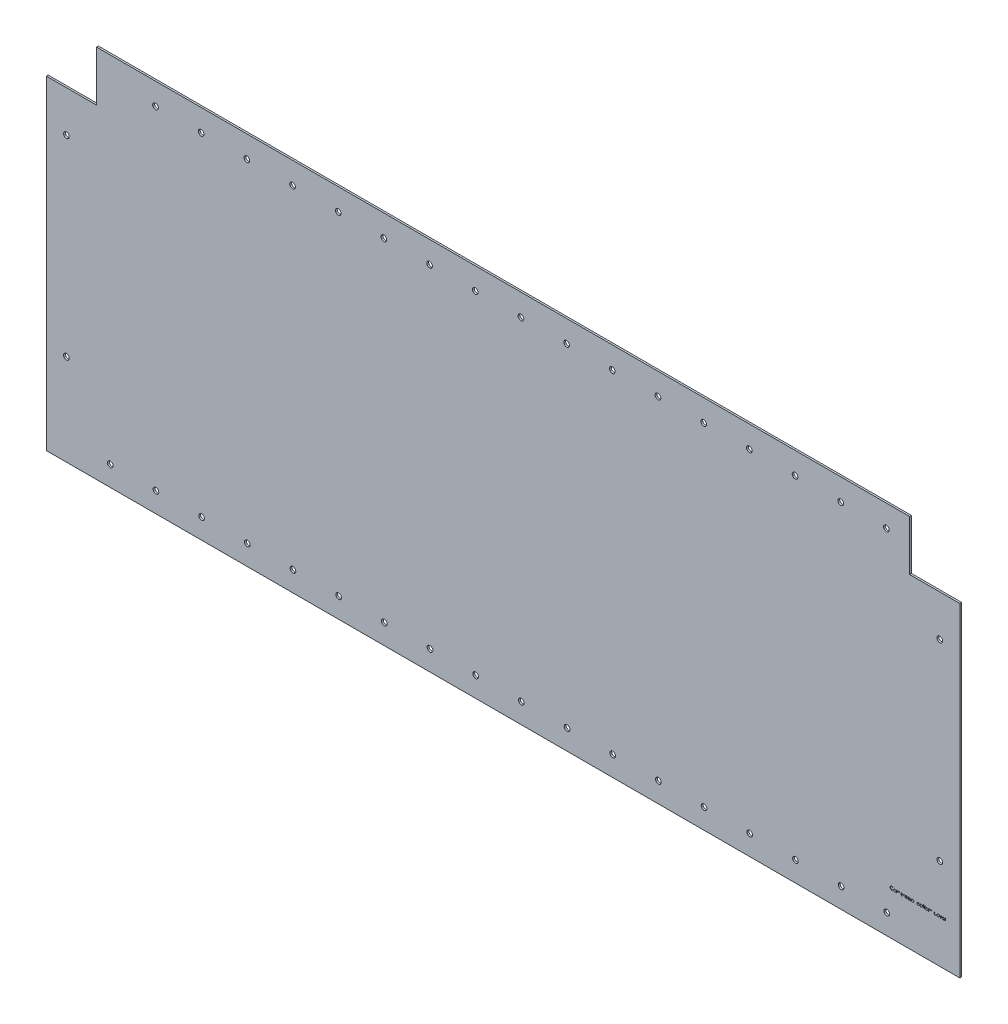
SolidWorks part; units mm, degrees
ref_plane "Front Plane" through (0, 0, 0) normal (0, 0, 1) x (1, 0, 0)
ref_plane "Top Plane" through (0, 0, 0) normal (0, 1, 0) x (1, 0, 0)
ref_plane "Right Plane" through (0, 0, 0) normal (1, 0, 0) x (0, 0, -1)
sketch "Sketch1" plane through (0, 0, 0) normal (0, 0, 1) x (1, 0, 0)
  line L0 (22, -100) -> (22, -380.8281) construction
  line L1 (0, 0) -> (1000, 0)
  line L2 (0, 0) -> (0, -410)
  line L3 (0, -410) -> (1000, -410)
  line L4 (1000, 0) -> (1000, -410)
  line L5 (22, -100) -> (940.6914, -100) construction
  line L6 (978, -100) -> (978, -347.1788) construction
  line L7 (22, -310) -> (989.4828, -310) construction
  circle A0 centre (22, -100) radius 3.1
  circle A1 centre (22, -310) radius 3.1
  circle A2 centre (978, -310) radius 3.1
  circle A3 centre (978, -100) radius 3.1
  dimension "D7" = 6.2
  dimension "D1" = 410
  dimension "D2" = 1000
  dimension "D3" = 22
  dimension "D4" = 100
  dimension "D5" = 100
  dimension "D6" = 22
extrude "Boss-Extrude1" add sketch "Sketch1" along normal blind 2
sketch "Sketch2" plane through (0, 0, 2) normal (0, 0, 1) x (1, 0, 0)
  line L0 (500, 0) -> (500, -410) construction
  line L1 (1000, 0) -> (945, 0)
  line L2 (1000, 0) -> (1000, -55)
  line L3 (1000, -55) -> (945, -55)
  line L4 (945, 0) -> (945, -55)
  line L5 (1000, 0) -> (0, 0) construction
  line L6 (0, -410) -> (1000, -410) construction
  line L7 (0, -55) -> (55, -55)
  line L8 (55, 0) -> (55, -55)
  line L9 (0, 0) -> (55, 0)
  line L10 (0, 0) -> (0, -55)
  dimension "D1" = 55
  dimension "D2" = 55
extrude "Cut-Extrude1" cut sketch "Sketch2" against normal blind 10
sketch "Sketch3" plane through (0, 0, 2) normal (0, 0, 1) x (1, 0, 0)
  line L0 (0, -388) -> (979.9055, -388) construction
  line L3 (0, -55) -> (0, -410) construction
  line L4 (0, -410) -> (1000, -410) construction
  circle A0 centre (70, -388) radius 3.1
  circle A1 centre (120, -388) radius 3.1
  circle A2 centre (170, -388) radius 3.1
  circle A3 centre (220, -388) radius 3.1
  circle A4 centre (270, -388) radius 3.1
  circle A5 centre (320, -388) radius 3.1
  circle A6 centre (370, -388) radius 3.1
  circle A7 centre (420, -388) radius 3.1
  circle A8 centre (470, -388) radius 3.1
  circle A9 centre (520, -388) radius 3.1
  circle A10 centre (570, -388) radius 3.1
  circle A11 centre (620, -388) radius 3.1
  circle A12 centre (670, -388) radius 3.1
  circle A13 centre (720, -388) radius 3.1
  circle A14 centre (770, -388) radius 3.1
  circle A15 centre (820, -388) radius 3.1
  circle A16 centre (870, -388) radius 3.1
  circle A17 centre (920, -388) radius 3.1
  dimension "D2" = 6.2
  dimension "D1" = 22
  dimension "D3" = 70
  dimension "D4" = 18
extrude "Cut-Extrude2" cut sketch "Sketch3" against normal through all
sketch "Sketch4" plane through (0, 0, 2) normal (0, 0, 1) x (1, 0, 0)
  line L0 (105, -24) -> (905.9107, -24) construction
  line L1 (945, 0) -> (55, 0) construction
  line L2 (55, -55) -> (55, 0) construction
  circle A0 centre (119.5493, -24) radius 3.1
  circle A1 centre (169.5493, -24) radius 3.1
  circle A2 centre (219.5493, -24) radius 3.1
  circle A3 centre (269.5493, -24) radius 3.1
  circle A4 centre (319.5493, -24) radius 3.1
  circle A5 centre (369.5493, -24) radius 3.1
  circle A6 centre (419.5493, -24) radius 3.1
  circle A7 centre (469.5493, -24) radius 3.1
  circle A8 centre (519.5493, -24) radius 3.1
  circle A9 centre (569.5493, -24) radius 3.1
  circle A10 centre (619.5493, -24) radius 3.1
  circle A11 centre (669.5493, -24) radius 3.1
  circle A12 centre (719.5493, -24) radius 3.1
  circle A13 centre (769.5493, -24) radius 3.1
  circle A14 centre (819.5493, -24) radius 3.1
  circle A15 centre (869.5493, -24) radius 3.1
  circle A16 centre (919.5493, -24) radius 3.1
  dimension "D3" = 6.2
  dimension "D1" = 24
  dimension "D2" = 50
  dimension "D4" = 17
extrude "Cut-Extrude3" cut sketch "Sketch4" against normal through all
sketch "Sketch5" plane through (0, 0, 2) normal (0, 0, 1) x (1, 0, 0)
  line L0 (923.3148, -363.8914) -> (994.2448, -363.8914) construction
  line L1 (926.9943, -361.0336) -> (926.7195, -361.244)
  line L2 (926.7195, -363.0388) -> (926.9943, -363.2471)
  line L3 (930.8084, -361.3337) -> (931.1225, -361.3337)
  line L4 (931.1225, -361.3337) -> (931.1225, -361.7782)
  line L5 (934.6225, -362.506) -> (934.6225, -363.8914)
  line L6 (934.6225, -363.8914) -> (934.3084, -363.8914)
  line L7 (934.3084, -363.8914) -> (934.3084, -362.5046)
  line L8 (932.8725, -362.8965) -> (932.8725, -363.8914)
  line L9 (932.8725, -363.8914) -> (932.5584, -363.8914)
  line L10 (932.5584, -363.8914) -> (932.5584, -362.5908)
  line L11 (931.1225, -362.8152) -> (931.1225, -363.8914)
  line L12 (931.1225, -363.8914) -> (930.8084, -363.8914)
  line L13 (930.8084, -363.8914) -> (930.8084, -361.3337)
  line L14 (935.3405, -361.3337) -> (935.6546, -361.3337)
  line L15 (935.6546, -361.3337) -> (935.6546, -361.807)
  line L16 (935.6546, -363.428) -> (935.6546, -364.8337)
  line L17 (935.6546, -364.8337) -> (935.3405, -364.8337)
  line L18 (935.3405, -364.8337) -> (935.3405, -361.3337)
  line L19 (938.5713, -361.3337) -> (938.8854, -361.3337)
  line L20 (938.8854, -361.3337) -> (938.8854, -361.7102)
  line L21 (939.7828, -361.3765) -> (939.6103, -361.6485)
  line L22 (938.8854, -363.0318) -> (938.8854, -363.8914)
  line L23 (938.8854, -363.8914) -> (938.5713, -363.8914)
  line L24 (938.5713, -363.8914) -> (938.5713, -361.3337)
  line L25 (942.1961, -363.0837) -> (942.4751, -363.2302)
  line L26 (942.6097, -362.6799) -> (940.3213, -362.6799)
  line L27 (940.3542, -362.3658) -> (942.2956, -362.3658)
  line L28 (944.4495, -361.6527) -> (944.2363, -361.8722)
  line L29 (943.0136, -363.5899) -> (943.2218, -363.3529)
  line L30 (946.3341, -361.6527) -> (946.1209, -361.8722)
  line L31 (944.8982, -363.5899) -> (945.1064, -363.3529)
  line L32 (950.1033, -361.3337) -> (950.4174, -361.3337)
  line L33 (950.4174, -361.3337) -> (950.4174, -361.7102)
  line L34 (951.3148, -361.3765) -> (951.1424, -361.6485)
  line L35 (950.4174, -363.0318) -> (950.4174, -363.8914)
  line L36 (950.4174, -363.8914) -> (950.1033, -363.8914)
  line L37 (950.1033, -363.8914) -> (950.1033, -361.3337)
  line L38 (952.9751, -363.8914) -> (952.9751, -360.3017)
  line L39 (952.9751, -360.3017) -> (953.2892, -360.3017)
  line L40 (953.2892, -360.3017) -> (953.2892, -361.7978)
  line L41 (953.2892, -363.4181) -> (953.2892, -363.8914)
  line L42 (953.2892, -363.8914) -> (952.9751, -363.8914)
  line L43 (959.7956, -360.3017) -> (960.1097, -360.3017)
  line L44 (960.1097, -360.3017) -> (960.1097, -361.3337)
  line L45 (960.1097, -361.3337) -> (960.5584, -361.3337)
  line L46 (960.5584, -361.3337) -> (960.5584, -361.6478)
  line L47 (960.5584, -361.6478) -> (960.1097, -361.6478)
  line L48 (960.1097, -361.6478) -> (960.1097, -363.8914)
  line L49 (960.1097, -363.8914) -> (959.7956, -363.8914)
  line L50 (959.7956, -363.8914) -> (959.7956, -361.6478)
  line L51 (959.7956, -361.6478) -> (959.3469, -361.6478)
  line L52 (959.3469, -361.6478) -> (959.3469, -361.3337)
  line L53 (959.3469, -361.3337) -> (959.7956, -361.3337)
  line L54 (959.7956, -361.3337) -> (959.7956, -360.3017)
  line L55 (961.411, -360.3017) -> (961.7251, -360.3017)
  line L56 (961.7251, -360.3017) -> (961.7251, -361.3337)
  line L57 (961.7251, -361.3337) -> (962.1738, -361.3337)
  line L58 (962.1738, -361.3337) -> (962.1738, -361.6478)
  line L59 (962.1738, -361.6478) -> (961.7251, -361.6478)
  line L60 (961.7251, -361.6478) -> (961.7251, -363.8914)
  line L61 (961.7251, -363.8914) -> (961.411, -363.8914)
  line L62 (961.411, -363.8914) -> (961.411, -361.6478)
  line L63 (961.411, -361.6478) -> (960.9623, -361.6478)
  line L64 (960.9623, -361.6478) -> (960.9623, -361.3337)
  line L65 (960.9623, -361.3337) -> (961.411, -361.3337)
  line L66 (961.411, -361.3337) -> (961.411, -360.3017)
  line L67 (965.8982, -361.3337) -> (966.2123, -361.3337)
  line L68 (966.2123, -361.3337) -> (966.2123, -361.7782)
  line L69 (969.7123, -362.506) -> (969.7123, -363.8914)
  line L70 (969.7123, -363.8914) -> (969.3982, -363.8914)
  line L71 (969.3982, -363.8914) -> (969.3982, -362.5046)
  line L72 (967.9623, -362.8965) -> (967.9623, -363.8914)
  line L73 (967.9623, -363.8914) -> (967.6482, -363.8914)
  line L74 (967.6482, -363.8914) -> (967.6482, -362.5908)
  line L75 (966.2123, -362.8152) -> (966.2123, -363.8914)
  line L76 (966.2123, -363.8914) -> (965.8982, -363.8914)
  line L77 (965.8982, -363.8914) -> (965.8982, -361.3337)
  line L78 (974.2892, -361.8883) -> (974.0263, -362.0517)
  line L79 (974.0263, -363.1734) -> (974.2892, -363.3459)
  line L80 (977.8341, -361.3337) -> (978.1741, -361.3337)
  line L81 (978.1741, -361.3337) -> (979.0232, -363.1959)
  line L82 (979.0232, -363.1959) -> (979.8722, -361.3337)
  line L83 (979.8722, -361.3337) -> (980.2123, -361.3337)
  line L84 (980.2123, -361.3337) -> (979.0456, -363.8914)
  line L85 (979.0456, -363.8914) -> (979.0007, -363.8914)
  line L86 (979.0007, -363.8914) -> (977.8341, -361.3337)
  line L87 (982.8499, -363.0837) -> (983.129, -363.2302)
  line L88 (983.2636, -362.6799) -> (980.9751, -362.6799)
  line L89 (981.0081, -362.3658) -> (982.9495, -362.3658)
  line L90 (983.802, -361.3337) -> (984.1161, -361.3337)
  line L91 (984.1161, -361.3337) -> (984.1161, -361.7102)
  line L92 (985.0136, -361.3765) -> (984.8411, -361.6485)
  line L93 (984.1161, -363.0318) -> (984.1161, -363.8914)
  line L94 (984.1161, -363.8914) -> (983.802, -363.8914)
  line L95 (983.802, -363.8914) -> (983.802, -361.3337)
  spline S0 degree 3 poles (926.7195, -361.244) (926.6812, -361.197) (926.6206, -361.1298) (926.533, -361.0479) (926.4651, -360.9907) (926.3933, -360.9393) (926.3194, -360.891) (926.2422, -360.8477) (926.1355, -360.7953) (925.9958, -360.7406) (925.7584, -360.6782) (925.5728, -360.66) (925.4477, -360.6606) knots 0 0 0 0 0.125475 0.187121 0.248294 0.309295 0.36985 0.430973 0.492456 0.616148 0.740844 1 1 1 1
  spline S1 degree 3 poles (925.4477, -360.6606) (925.3778, -360.6597) (925.2738, -360.6672) (925.1374, -360.6874) (925.0377, -360.7095) (924.9401, -360.7375) (924.844, -360.7709) (924.7508, -360.8122) (924.6592, -360.8579) (924.5714, -360.9096) (924.4883, -360.9659) (924.4103, -361.0263) (924.3372, -361.0909) (924.2691, -361.1595) (924.2063, -361.2329) (924.1491, -361.3108) (924.0964, -361.3921) (924.0492, -361.4766) (924.0096, -361.5647) (923.9746, -361.6548) (923.9469, -361.7479) (923.925, -361.8435) (923.9045, -361.9757) (923.8973, -362.0767) (923.8982, -362.1449) knots 0 0 0 0 0.087502 0.130463 0.172752 0.215403 0.25765 0.300153 0.343121 0.385925 0.427686 0.468818 0.509492 0.549883 0.58998 0.630405 0.670869 0.711384 0.751627 0.791776 0.832459 0.873319 0.914543 1 1 1 1
  spline S2 degree 3 poles (923.8982, -362.1449) (923.8977, -362.2465) (923.9119, -362.3966) (923.9575, -362.5895) (924.0077, -362.7249) (924.0696, -362.8548) (924.1478, -362.977) (924.2385, -363.0934) (924.3427, -363.2013) (924.4571, -363.2998) (924.5799, -363.3865) (924.7107, -363.4589) (924.8481, -363.519) (924.9931, -363.5652) (925.1998, -363.6097) (925.3604, -363.623) (925.4694, -363.6222) knots 0 0 0 0 0.12629 0.186726 0.246146 0.305576 0.365429 0.426326 0.48884 0.551725 0.613919 0.675484 0.737334 0.800229 0.864502 1 1 1 1
  spline S3 degree 3 poles (925.4694, -363.6222) (925.5896, -363.6222) (925.7681, -363.6053) (925.996, -363.5433) (926.1573, -363.4795) (926.3106, -363.3963) (926.5082, -363.26) (926.6388, -363.1317) (926.7195, -363.0388) knots 0 0 0 0 0.252949 0.374755 0.49594 0.617181 0.740909 1 1 1 1
  spline S4 degree 3 poles (926.9943, -363.2471) (926.951, -363.3046) (926.8822, -363.3873) (926.7813, -363.4883) (926.7017, -363.5585) (926.6186, -363.6246) (926.5305, -363.6849) (926.4386, -363.7402) (926.3433, -363.7908) (926.2445, -363.8357) (926.1425, -363.8742) (926.0377, -363.9073) (925.93, -363.9346) (925.8193, -363.9558) (925.6665, -363.9751) (925.55, -363.9817) (925.4715, -363.9811) knots 0 0 0 0 0.123053 0.183475 0.243727 0.304279 0.364863 0.425946 0.487391 0.54922 0.611144 0.673529 0.736961 0.800785 0.866013 1 1 1 1
  spline S5 degree 3 poles (925.4715, -363.9811) (925.397, -363.9821) (925.2869, -363.9761) (925.1425, -363.9605) (925.0388, -363.9433) (924.9376, -363.9229) (924.8401, -363.8957) (924.7451, -363.8651) (924.6531, -363.8292) (924.5641, -363.7887) (924.4782, -363.7429) (924.3956, -363.6922) (924.3154, -363.6378) (924.2388, -363.5778) (924.1399, -363.4911) (924.071, -363.4197) (924.0279, -363.3691) knots 0 0 0 0 0.13775 0.203917 0.26878 0.332414 0.394754 0.45618 0.516996 0.577396 0.637198 0.696999 0.756756 0.816554 0.876948 1 1 1 1
  spline S6 degree 3 poles (924.0279, -363.3691) (923.9554, -363.2843) (923.8579, -363.1485) (923.7548, -362.9522) (923.6923, -362.7988) (923.6436, -362.6388) (923.5977, -362.4133) (923.5837, -362.2389) (923.5841, -362.1211) knots 0 0 0 0 0.247156 0.36878 0.490734 0.613614 0.738958 1 1 1 1
  spline S7 degree 3 poles (923.5841, -362.1211) (923.584, -361.9973) (923.5997, -361.8138) (923.6566, -361.5783) (923.7159, -361.4121) (923.7912, -361.253) (923.8842, -361.1021) (923.9939, -360.9586) (924.1194, -360.8246) (924.2569, -360.7021) (924.4042, -360.5943) (924.561, -360.5046) (924.7255, -360.4295) (924.899, -360.372) (925.1456, -360.317) (925.3375, -360.3019) (925.4673, -360.3017) knots 0 0 0 0 0.127014 0.187955 0.248014 0.307748 0.368235 0.42947 0.492743 0.556258 0.618217 0.679655 0.741246 0.803415 0.866815 1 1 1 1
  spline S8 degree 3 poles (925.4673, -360.3017) (925.5469, -360.3015) (925.665, -360.3069) (925.8195, -360.3279) (925.9311, -360.349) (926.0402, -360.3752) (926.146, -360.4094) (926.2491, -360.4484) (926.3489, -360.4934) (926.4448, -360.5438) (926.5369, -360.5993) (926.6243, -360.6595) (926.7078, -360.7242) (926.7859, -360.7946) (926.8862, -360.8938) (926.9521, -360.9769) (926.9943, -361.0336) knots 0 0 0 0 0.135683 0.201215 0.265682 0.329267 0.392395 0.45507 0.517127 0.57879 0.63974 0.700192 0.759806 0.819628 0.879355 1 1 1 1
  spline S9 degree 3 poles (928.8579, -361.2888) (928.952, -361.2879) (929.0912, -361.3014) (929.2694, -361.3461) (929.3952, -361.3913) (929.5135, -361.452) (929.6659, -361.5495) (929.7675, -361.6423) (929.8297, -361.7102) knots 0 0 0 0 0.258332 0.382134 0.503804 0.624693 0.746871 1 1 1 1
  spline S10 degree 3 poles (929.8297, -361.7102) (929.8867, -361.7725) (929.9631, -361.8725) (930.0453, -362.0168) (930.0944, -362.1291) (930.1331, -362.2454) (930.1703, -362.4084) (930.1798, -362.5346) (930.1802, -362.6196) knots 0 0 0 0 0.253834 0.376506 0.498534 0.621368 0.744565 1 1 1 1
  spline S11 degree 3 poles (930.1802, -362.6196) (930.1807, -362.7051) (930.169, -362.8323) (930.1304, -362.9966) (930.0896, -363.1145) (930.0372, -363.2284) (929.9734, -363.3378) (929.8975, -363.4429) (929.8115, -363.5429) (929.7164, -363.6351) (929.6133, -363.7154) (929.5042, -363.7843) (929.3875, -363.8397) (929.2644, -363.8834) (929.0884, -363.9252) (928.9509, -363.9359) (928.8579, -363.9363) knots 0 0 0 0 0.123337 0.183265 0.243172 0.302898 0.363774 0.425605 0.489659 0.553785 0.616222 0.677854 0.739517 0.802097 0.865866 1 1 1 1
  spline S12 degree 3 poles (928.8579, -363.9363) (928.7645, -363.9358) (928.6265, -363.9254) (928.45, -363.8834) (928.3267, -363.8396) (928.2096, -363.7843) (928.0998, -363.7156) (927.9966, -363.6351) (927.9015, -363.543) (927.8155, -363.4429) (927.7397, -363.3378) (927.6758, -363.2284) (927.6234, -363.1145) (927.5826, -362.9966) (927.544, -362.8323) (927.5323, -362.7051) (927.5328, -362.6196) knots 0 0 0 0 0.134635 0.198324 0.260825 0.322714 0.384555 0.446913 0.510958 0.574931 0.636685 0.697483 0.757134 0.816966 0.876818 1 1 1 1
  spline S13 degree 3 poles (927.5328, -362.6196) (927.5333, -362.5349) (927.5428, -362.4089) (927.5799, -362.2464) (927.6185, -362.1304) (927.6681, -362.0187) (927.7492, -361.8739) (927.8269, -361.7748) (927.8834, -361.7123) knots 0 0 0 0 0.255238 0.378679 0.501088 0.622714 0.746241 1 1 1 1
  spline S14 degree 3 poles (927.8834, -361.7123) (927.945, -361.6435) (928.0475, -361.5516) (928.1995, -361.4521) (928.3192, -361.3926) (928.4449, -361.3458) (928.6237, -361.3015) (928.7633, -361.288) (928.8579, -361.2888) knots 0 0 0 0 0.252713 0.374819 0.496436 0.617911 0.741288 1 1 1 1
  spline S15 degree 3 poles (928.8565, -361.6029) (928.7895, -361.6031) (928.69, -361.6122) (928.562, -361.6433) (928.4706, -361.6758) (928.3829, -361.7179) (928.299, -361.7696) (928.2186, -361.8303) (928.1432, -361.8997) (928.074, -361.9756) (928.0136, -362.0565) (927.9621, -362.141) (927.9193, -362.2292) (927.8874, -362.3221) (927.856, -362.4523) (927.8471, -362.5535) (927.8469, -362.6217) knots 0 0 0 0 0.126044 0.187165 0.247399 0.30838 0.36978 0.432584 0.497641 0.562401 0.625557 0.687332 0.748313 0.809791 0.871768 1 1 1 1
  spline S16 degree 3 poles (927.8469, -362.6217) (927.8471, -362.7104) (927.8627, -362.8437) (927.9211, -363.0116) (927.9796, -363.1313) (928.053, -363.2419) (928.1395, -363.3406) (928.2381, -363.4258) (928.3478, -363.4965) (928.4661, -363.5526) (928.6345, -363.6064) (928.7672, -363.6232) (928.8565, -363.6222) knots 0 0 0 0 0.168179 0.251488 0.335841 0.419834 0.502345 0.583649 0.665931 0.748717 0.831047 1 1 1 1
  spline S17 degree 3 poles (928.8565, -363.6222) (928.9458, -363.6231) (929.0784, -363.6067) (929.2464, -363.5524) (929.3646, -363.4965) (929.4742, -363.4255) (929.5735, -363.3411) (929.6593, -363.2417) (929.7326, -363.1311) (929.7921, -363.0118) (929.8502, -362.8436) (929.866, -362.7104) (929.8661, -362.6217) knots 0 0 0 0 0.168983 0.250908 0.333708 0.416005 0.49766 0.579893 0.663902 0.748466 0.831791 1 1 1 1
  spline S18 degree 3 poles (929.8661, -362.6217) (929.8659, -362.5535) (929.857, -362.4523) (929.8256, -362.3221) (929.7937, -362.2293) (929.751, -362.1407) (929.6986, -362.0567) (929.6384, -361.9753) (929.5684, -361.9) (929.4931, -361.8303) (929.4126, -361.7696) (929.3288, -361.7182) (929.2414, -361.6755) (929.15, -361.6436) (929.0224, -361.6119) (928.9232, -361.6033) (928.8565, -361.6029) knots 0 0 0 0 0.128274 0.19027 0.251768 0.312769 0.374793 0.43797 0.503047 0.568125 0.63095 0.692369 0.752973 0.813641 0.874355 1 1 1 1
  spline S19 degree 3 poles (931.1225, -361.7782) (931.1752, -361.7028) (931.2816, -361.5699) (931.4116, -361.4598) (931.4773, -361.4185) knots 0 0 0 0 0.543395 1 1 1 1
  spline S20 degree 3 poles (931.4773, -361.4185) (931.5589, -361.3764) (931.7307, -361.3097) (931.9138, -361.2895) (932.0046, -361.2888) knots 0 0 0 0 0.503035 1 1 1 1
  spline S21 degree 3 poles (932.0046, -361.2888) (932.0656, -361.2896) (932.1572, -361.2974) (932.275, -361.3287) (932.3596, -361.3611) (932.4394, -361.4003) (932.5124, -361.4464) (932.5781, -361.4981) (932.6362, -361.5578) (932.6885, -361.6271) (932.7562, -361.7409) (932.795, -361.8379) (932.8186, -361.9065) knots 0 0 0 0 0.166532 0.248836 0.331246 0.412957 0.490494 0.566156 0.639987 0.716765 0.802144 1 1 1 1
  spline S22 degree 3 poles (932.8186, -361.9065) (932.8447, -361.8574) (932.8877, -361.787) (932.952, -361.6999) (933.0021, -361.6399) (933.0545, -361.5846) (933.1095, -361.5338) (933.1669, -361.4873) (933.2467, -361.4329) (933.3505, -361.3753) (933.5251, -361.3082) (933.6643, -361.2886) (933.7567, -361.2888) knots 0 0 0 0 0.141226 0.209116 0.27484 0.339483 0.402476 0.464942 0.526833 0.647415 0.765562 1 1 1 1
  spline S23 degree 3 poles (933.7567, -361.2888) (933.8403, -361.2895) (933.9653, -361.3032) (934.1196, -361.3612) (934.2251, -361.4194) (934.3202, -361.4926) (934.4029, -361.5796) (934.4727, -361.68) (934.5183, -361.7744) (934.5492, -361.8577) (934.5683, -361.9287) (934.5851, -362.0069) (934.5991, -362.0922) (934.6093, -362.1852) (934.6198, -362.3237) (934.6229, -362.4316) (934.6225, -362.506) knots 0 0 0 0 0.147965 0.218797 0.28947 0.359724 0.429708 0.500497 0.574429 0.613947 0.657155 0.703973 0.754939 0.809707 0.868833 1 1 1 1
  spline S24 degree 3 poles (934.3084, -362.5046) (934.3085, -362.4417) (934.3075, -362.3514) (934.3004, -362.2365) (934.2945, -362.1623) (934.2863, -362.096) (934.2756, -362.0378) (934.2643, -361.9872) (934.2456, -361.9312) (934.2157, -361.8693) (934.17, -361.8026) (934.1126, -361.7445) (934.0462, -361.6941) (933.9707, -361.6531) (933.8568, -361.6129) (933.7645, -361.6025) (933.702, -361.6029) knots 0 0 0 0 0.150563 0.216151 0.27568 0.328707 0.375904 0.417302 0.452693 0.517265 0.581217 0.645322 0.712024 0.78013 0.850218 1 1 1 1
  spline S25 degree 3 poles (933.702, -361.6029) (933.6234, -361.6016) (933.5064, -361.6209) (933.3595, -361.6789) (933.2573, -361.7412) (933.1632, -361.8161) (933.0823, -361.905) (933.0155, -362.0056) (932.9702, -362.0988) (932.9417, -362.1824) (932.9228, -362.2555) (932.9081, -362.3386) (932.8943, -362.4311) (932.8853, -362.5337) (932.874, -362.6897) (932.873, -362.8119) (932.8725, -362.8965) knots 0 0 0 0 0.134707 0.201865 0.270788 0.340024 0.408083 0.476813 0.547346 0.58564 0.628865 0.677153 0.730803 0.789807 0.854325 1 1 1 1
  spline S26 degree 3 poles (932.5584, -362.5908) (932.5585, -362.5202) (932.5576, -362.4189) (932.5504, -362.2902) (932.5446, -362.2074) (932.5361, -362.134) (932.5265, -362.0696) (932.5151, -362.0144) (932.4964, -361.9538) (932.4676, -361.8871) (932.4215, -361.8159) (932.3638, -361.7537) (932.2963, -361.7005) (932.2203, -361.6566) (932.1059, -361.6133) (932.0125, -361.6035) (931.9499, -361.6029) knots 0 0 0 0 0.158779 0.227738 0.289946 0.345499 0.393896 0.436374 0.472122 0.536384 0.599078 0.661948 0.726311 0.791771 0.858647 1 1 1 1
  spline S27 degree 3 poles (931.9499, -361.6029) (931.8741, -361.6023) (931.7601, -361.6205) (931.6173, -361.678) (931.5153, -361.7376) (931.4217, -361.8115) (931.3397, -361.8984) (931.2707, -361.9973) (931.225, -362.0895) (931.1955, -362.171) (931.1759, -362.2404) (931.1591, -362.3174) (931.1465, -362.4023) (931.1345, -362.4945) (931.1263, -362.633) (931.1215, -362.7408) (931.1225, -362.8152) knots 0 0 0 0 0.136871 0.206114 0.277538 0.349772 0.421251 0.492911 0.567027 0.606614 0.649704 0.697303 0.749086 0.804881 0.865485 1 1 1 1
  spline S28 degree 3 poles (935.6546, -361.807) (935.7168, -361.7217) (935.8212, -361.6057) (935.9825, -361.4815) (936.1096, -361.4101) (936.244, -361.3564) (936.4352, -361.3022) (936.5863, -361.2892) (936.688, -361.2888) knots 0 0 0 0 0.263045 0.386061 0.505771 0.625178 0.746148 1 1 1 1
  spline S29 degree 3 poles (936.688, -361.2888) (936.7777, -361.2897) (936.911, -361.2997) (937.0824, -361.3405) (937.204, -361.3838) (937.3212, -361.4375) (937.4324, -361.5052) (937.5394, -361.5836) (937.6393, -361.6738) (937.7316, -361.7715) (937.8114, -361.8765) (937.8803, -361.9855) (937.936, -362.1) (937.9796, -362.2194) (938.0215, -362.3871) (938.0323, -362.5177) (938.0328, -362.6055) knots 0 0 0 0 0.128636 0.190653 0.252125 0.313446 0.375227 0.438498 0.503285 0.56801 0.630879 0.692154 0.752552 0.813191 0.873985 1 1 1 1
  spline S30 degree 3 poles (938.0328, -362.6055) (938.0326, -362.695) (938.0211, -362.8277) (937.9804, -362.9985) (937.9374, -363.1197) (937.8818, -363.2357) (937.814, -363.3463) (937.7342, -363.4515) (937.6429, -363.5499) (937.5438, -363.6405) (937.4379, -363.7197) (937.3269, -363.7862) (937.2112, -363.8418) (937.0899, -363.8837) (936.9196, -363.9246) (936.7871, -363.9359) (936.6979, -363.9363) knots 0 0 0 0 0.128034 0.189574 0.25058 0.311733 0.37325 0.435763 0.500346 0.564949 0.627528 0.689157 0.749865 0.81076 0.8723 1 1 1 1
  spline S31 degree 3 poles (936.6979, -363.9363) (936.5974, -363.9374) (936.4489, -363.9203) (936.2586, -363.8677) (936.1244, -363.8111) (935.9962, -363.7388) (935.8312, -363.6193) (935.7221, -363.5081) (935.6546, -363.428) knots 0 0 0 0 0.250548 0.37123 0.492116 0.613401 0.737997 1 1 1 1
  spline S32 degree 3 poles (936.6852, -361.6029) (936.6151, -361.6019) (936.5117, -361.612) (936.378, -361.6416) (936.2839, -361.6745) (936.1937, -361.7149) (936.108, -361.7653) (936.0269, -361.825) (935.9507, -361.8927) (935.8818, -361.9672) (935.8209, -362.0468) (935.7697, -362.1313) (935.7272, -362.22) (935.6949, -362.3134) (935.6636, -362.4456) (935.6548, -362.5486) (935.6546, -362.6182) knots 0 0 0 0 0.130024 0.192374 0.253884 0.314896 0.375806 0.438242 0.501591 0.564881 0.626533 0.687516 0.748106 0.808796 0.870822 1 1 1 1
  spline S33 degree 3 poles (935.6546, -362.6182) (935.6548, -362.7089) (935.6699, -362.844) (935.7259, -363.0139) (935.7844, -363.1313) (935.8584, -363.2393) (935.9474, -363.336) (936.0509, -363.4208) (936.167, -363.4922) (936.2914, -363.5501) (936.4645, -363.6059) (936.6, -363.622) (936.6901, -363.6222) knots 0 0 0 0 0.169344 0.251061 0.332326 0.413189 0.494299 0.576654 0.661785 0.747765 0.831967 1 1 1 1
  spline S34 degree 3 poles (936.6901, -363.6222) (936.7786, -363.6227) (936.9108, -363.6048) (937.0797, -363.5499) (937.1999, -363.4904) (937.3127, -363.4174) (937.4146, -363.3298) (937.5036, -363.2283) (937.5795, -363.1153) (937.6406, -362.9942) (937.7018, -362.8277) (937.7177, -362.6959) (937.7187, -362.609) knots 0 0 0 0 0.165574 0.248159 0.332033 0.416257 0.499525 0.583039 0.668596 0.754035 0.83692 1 1 1 1
  spline S35 degree 3 poles (937.7187, -362.609) (937.7199, -362.5215) (937.7003, -362.3906) (937.6428, -362.2232) (937.5804, -362.1036) (937.5061, -361.9909) (937.4164, -361.8913) (937.3158, -361.8042) (937.2031, -361.7321) (937.0821, -361.6749) (936.9111, -361.6183) (936.7757, -361.6033) (936.6852, -361.6029) knots 0 0 0 0 0.163349 0.245826 0.330367 0.415198 0.497941 0.580476 0.66374 0.747513 0.830399 1 1 1 1
  spline S36 degree 3 poles (938.8854, -361.7102) (938.9284, -361.6425) (938.9963, -361.5487) (939.1021, -361.446) (939.1798, -361.3875) (939.2601, -361.3437) (939.3677, -361.3011) (939.4533, -361.2892) (939.5094, -361.2888) knots 0 0 0 0 0.306112 0.438367 0.560541 0.675317 0.786114 1 1 1 1
  spline S37 degree 3 poles (939.5094, -361.2888) (939.5543, -361.2892) (939.6508, -361.3061) (939.7385, -361.3496) (939.7828, -361.3765) knots 0 0 0 0 0.463523 1 1 1 1
  spline S38 degree 3 poles (939.6103, -361.6485) (939.5817, -361.6358) (939.5302, -361.6126) (939.4744, -361.6033) (939.4498, -361.6029) knots 0 0 0 0 0.56023 1 1 1 1
  spline S39 degree 3 poles (939.4498, -361.6029) (939.3982, -361.6029) (939.3194, -361.6217) (939.2244, -361.6786) (939.1662, -361.7268) (939.1212, -361.7733) (939.0891, -361.814) (939.0596, -361.8596) (939.0314, -361.9093) (939.0057, -361.964) (938.9729, -362.0451) (938.9534, -362.1095) (938.9415, -362.154) knots 0 0 0 0 0.191338 0.295191 0.410312 0.47193 0.536425 0.603119 0.674118 0.749332 0.828283 1 1 1 1
  spline S40 degree 3 poles (938.9415, -362.154) (938.9297, -362.1987) (938.9182, -362.2738) (938.906, -362.3836) (938.8989, -362.4865) (938.8923, -362.6031) (938.887, -362.7864) (938.8848, -362.9308) (938.8854, -363.0318) knots 0 0 0 0 0.156938 0.2586 0.375891 0.508166 0.656238 1 1 1 1
  spline S41 degree 3 poles (942.4751, -363.2302) (942.4336, -363.3079) (942.3641, -363.4169) (942.2572, -363.5467) (942.1721, -363.6284) (942.0824, -363.6997) (941.9877, -363.762) (941.8874, -363.8151) (941.7816, -363.8599) (941.6693, -363.8943) (941.5069, -363.9276) (941.38, -363.9363) (941.2937, -363.9363) knots 0 0 0 0 0.181661 0.265874 0.346355 0.4246 0.501903 0.579992 0.658443 0.738672 0.821894 1 1 1 1
  spline S42 degree 3 poles (941.2937, -363.9363) (941.1979, -363.9362) (941.057, -363.9252) (940.8778, -363.8821) (940.7546, -363.8382) (940.6398, -363.7807) (940.5333, -363.7108) (940.4345, -363.6286) (940.3465, -363.5336) (940.2672, -363.4319) (940.1973, -363.326) (940.1389, -363.216) (940.0913, -363.1027) (940.0529, -362.9869) (940.0168, -362.8264) (940.0081, -362.7026) (940.0072, -362.6196) knots 0 0 0 0 0.139629 0.204797 0.268135 0.329814 0.391301 0.453434 0.516552 0.579631 0.641119 0.701294 0.76081 0.819932 0.87892 1 1 1 1
  spline S43 degree 3 poles (940.0072, -362.6196) (940.0081, -362.5418) (940.0154, -362.4256) (940.047, -362.2751) (940.0792, -362.1662) (940.1207, -362.0607) (940.1889, -361.9232) (940.2541, -361.8271) (940.3016, -361.7656) knots 0 0 0 0 0.253768 0.377428 0.500551 0.623296 0.746578 1 1 1 1
  spline S44 degree 3 poles (940.3016, -361.7656) (940.3622, -361.6899) (940.461, -361.584) (940.6156, -361.4732) (940.7372, -361.4052) (940.8675, -361.3536) (941.0541, -361.3011) (941.202, -361.29) (941.3014, -361.2888) knots 0 0 0 0 0.253589 0.374643 0.49534 0.616325 0.739759 1 1 1 1
  spline S45 degree 3 poles (941.3014, -361.2888) (941.4043, -361.2884) (941.5562, -361.3033) (941.7488, -361.3566) (941.8826, -361.4117) (942.0083, -361.4829) (942.1665, -361.6019) (942.27, -361.7116) (942.3314, -361.7922) knots 0 0 0 0 0.259033 0.38188 0.502258 0.622752 0.744743 1 1 1 1
  spline S46 degree 3 poles (942.3314, -361.7922) (942.3773, -361.8511) (942.4372, -361.9468) (942.5008, -362.0836) (942.5392, -362.1924) (942.5702, -362.3063) (942.6008, -362.4686) (942.6081, -362.5946) (942.6097, -362.6799) knots 0 0 0 0 0.236255 0.356174 0.47725 0.60154 0.729618 1 1 1 1
  spline S47 degree 3 poles (940.3213, -362.6799) (940.323, -362.7461) (940.3319, -362.844) (940.3622, -362.9692) (940.3935, -363.0563) (940.4313, -363.1392) (940.4777, -363.2173) (940.5331, -363.2904) (940.5948, -363.359) (940.6635, -363.42) (940.7358, -363.4747) (940.8127, -363.5205) (940.8936, -363.5577) (940.9783, -363.5867) (941.0983, -363.6138) (941.1914, -363.6225) (941.2545, -363.6222) knots 0 0 0 0 0.134476 0.198391 0.260753 0.321829 0.383037 0.444653 0.507398 0.569825 0.630778 0.690929 0.750945 0.811049 0.872331 1 1 1 1
  spline S48 degree 3 poles (941.2545, -363.6222) (941.3166, -363.6225) (941.4099, -363.6151) (941.5318, -363.5896) (941.6211, -363.5638) (941.7066, -363.5322) (941.7859, -363.4941) (941.8587, -363.4519) (941.9269, -363.4037) (941.9929, -363.3447) (942.0864, -363.2399) (942.1535, -363.1503) (942.1961, -363.0837) knots 0 0 0 0 0.163879 0.245659 0.327726 0.40861 0.485749 0.559169 0.630268 0.705306 0.792065 1 1 1 1
  spline S49 degree 3 poles (942.2956, -362.3658) (942.2757, -362.285) (942.2361, -362.1711) (942.1637, -362.0342) (942.1021, -361.9486) (942.0322, -361.8726) (941.9516, -361.8062) (941.8612, -361.7468) (941.7614, -361.6966) (941.6558, -361.654) (941.508, -361.6154) (941.394, -361.6018) (941.3176, -361.6029) knots 0 0 0 0 0.185231 0.267501 0.3444 0.419595 0.496891 0.576638 0.660268 0.745387 0.83004 1 1 1 1
  spline S50 degree 3 poles (941.3176, -361.6029) (941.2556, -361.6028) (941.1636, -361.6095) (941.0453, -361.6352) (940.9605, -361.6611) (940.8799, -361.6958) (940.7749, -361.7502) (940.704, -361.8044) (940.6585, -361.8427) knots 0 0 0 0 0.259141 0.384162 0.505992 0.629098 0.750669 1 1 1 1
  spline S51 degree 3 poles (940.6585, -361.8427) (940.6236, -361.8721) (940.5764, -361.923) (940.5197, -361.9978) (940.4803, -362.0608) (940.4443, -362.1294) (940.398, -362.23) (940.3706, -362.3104) (940.3542, -362.3658) knots 0 0 0 0 0.22258 0.3385 0.458709 0.585535 0.717518 1 1 1 1
  spline S52 degree 3 poles (944.2363, -361.8722) (944.2015, -361.8306) (944.148, -361.7727) (944.0702, -361.7087) (944.0152, -361.6697) (943.9597, -361.6403) (943.8877, -361.6121) (943.8314, -361.603) (943.7946, -361.6029) knots 0 0 0 0 0.305036 0.441309 0.565963 0.683525 0.793334 1 1 1 1
  spline S53 degree 3 poles (943.7946, -361.6029) (943.751, -361.602) (943.6859, -361.6161) (943.6085, -361.6597) (943.5584, -361.7056) (943.5159, -361.7584) (943.4742, -361.8372) (943.4624, -361.9032) (943.4623, -361.9472) knots 0 0 0 0 0.245901 0.369166 0.498511 0.628504 0.751028 1 1 1 1
  spline S54 degree 3 poles (943.4623, -361.9472) (943.4624, -361.9876) (943.478, -362.0717) (943.5225, -362.1447) (943.5492, -362.1793) knots 0 0 0 0 0.479403 1 1 1 1
  spline S55 degree 3 poles (943.5492, -362.1793) (943.5652, -362.201) (943.5964, -362.2305) (943.642, -362.2707) (943.6853, -362.3027) (943.734, -362.3363) (943.8109, -362.3837) (943.8711, -362.4203) (943.9145, -362.4429) knots 0 0 0 0 0.17756 0.283982 0.402217 0.533568 0.676121 1 1 1 1
  spline S56 degree 3 poles (943.9145, -362.4429) (943.9672, -362.472) (944.0431, -362.5159) (944.1368, -362.5787) (944.1982, -362.6234) (944.2521, -362.6685) (944.3138, -362.7247) (944.353, -362.7706) (944.3751, -362.8019) knots 0 0 0 0 0.307115 0.446213 0.574876 0.694152 0.804581 1 1 1 1
  spline S57 degree 3 poles (944.3751, -362.8019) (944.4132, -362.8594) (944.4773, -362.986) (944.4933, -363.127) (944.4943, -363.1973) knots 0 0 0 0 0.495235 1 1 1 1
  spline S58 degree 3 poles (944.4943, -363.1973) (944.4939, -363.247) (944.4884, -363.3211) (944.4654, -363.4158) (944.4423, -363.4835) (944.4111, -363.5475) (944.3746, -363.6093) (944.3307, -363.6677) (944.2806, -363.7225) (944.2257, -363.7726) (944.1672, -363.8166) (944.105, -363.8532) (944.0395, -363.8835) (943.9705, -363.9075) (943.8725, -363.9302) (943.7962, -363.9359) (943.7448, -363.9363) knots 0 0 0 0 0.127199 0.188597 0.24864 0.309525 0.370037 0.431889 0.495704 0.559519 0.621372 0.682397 0.743568 0.805498 0.86864 1 1 1 1
  spline S59 degree 3 poles (943.7448, -363.9363) (943.6746, -363.9368) (943.5694, -363.9247) (943.4338, -363.886) (943.3354, -363.8463) (943.2424, -363.7961) (943.1292, -363.7165) (943.0558, -363.6435) (943.0136, -363.5899) knots 0 0 0 0 0.251724 0.377219 0.504694 0.631458 0.755401 1 1 1 1
  spline S60 degree 3 poles (943.2218, -363.3529) (943.2594, -363.3948) (943.3177, -363.4535) (943.4036, -363.517) (943.4664, -363.5557) (943.5306, -363.5854) (943.6171, -363.6133) (943.6843, -363.6224) (943.7287, -363.6222) knots 0 0 0 0 0.285904 0.417172 0.540501 0.659238 0.775006 1 1 1 1
  spline S61 degree 3 poles (943.7287, -363.6222) (943.7879, -363.6227) (943.8757, -363.6074) (943.9814, -363.5556) (944.0495, -363.5016) (944.1073, -363.4386) (944.1634, -363.3443) (944.1806, -363.2638) (944.1802, -363.2106) knots 0 0 0 0 0.261896 0.387836 0.517686 0.644509 0.764718 1 1 1 1
  spline S62 degree 3 poles (944.1802, -363.2106) (944.1801, -363.1666) (944.1661, -363.0783) (944.1219, -363.0006) (944.094, -362.9666) knots 0 0 0 0 0.500453 1 1 1 1
  spline S63 degree 3 poles (944.094, -362.9666) (944.0771, -362.9464) (944.0459, -362.9169) (943.998, -362.8789) (943.9529, -362.8465) (943.9009, -362.8129) (943.8183, -362.7643) (943.7526, -362.7275) (943.7063, -362.703) knots 0 0 0 0 0.167462 0.27227 0.389551 0.520801 0.666263 1 1 1 1
  spline S64 degree 3 poles (943.7063, -362.703) (943.6557, -362.675) (943.5827, -362.6333) (943.4936, -362.5717) (943.4345, -362.5288) (943.3824, -362.4853) (943.3245, -362.429) (943.2862, -362.3849) (943.2653, -362.3538) knots 0 0 0 0 0.30595 0.443775 0.572824 0.692154 0.802296 1 1 1 1
  spline S65 degree 3 poles (943.2653, -362.3538) (943.226, -362.2974) (943.1676, -362.1695) (943.1469, -362.0305) (943.1482, -361.9598) knots 0 0 0 0 0.492591 1 1 1 1
  spline S66 degree 3 poles (943.1482, -361.9598) (943.1485, -361.9137) (943.1526, -361.845) (943.1733, -361.7575) (943.1923, -361.6953) (943.2188, -361.6368) (943.2505, -361.5812) (943.2877, -361.5284) (943.3305, -361.4794) (943.3776, -361.4349) (943.4285, -361.3961) (943.4821, -361.363) (943.5385, -361.3352) (943.5983, -361.3143) (943.6835, -361.2945) (943.7497, -361.2883) (943.7946, -361.2888) knots 0 0 0 0 0.133044 0.196507 0.258613 0.319728 0.380873 0.442636 0.505079 0.567881 0.628814 0.68891 0.748765 0.809386 0.870884 1 1 1 1
  spline S67 degree 3 poles (943.7946, -361.2888) (943.8495, -361.2889) (943.9334, -361.3006) (944.0413, -361.339) (944.1236, -361.3792) (944.2054, -361.4313) (944.3189, -361.5182) (944.3989, -361.5954) (944.4495, -361.6527) knots 0 0 0 0 0.213412 0.326127 0.444452 0.569061 0.702712 1 1 1 1
  spline S68 degree 3 poles (946.1209, -361.8722) (946.0861, -361.8306) (946.0327, -361.7727) (945.9548, -361.7087) (945.8998, -361.6697) (945.8443, -361.6403) (945.7723, -361.6121) (945.716, -361.603) (945.6792, -361.6029) knots 0 0 0 0 0.305036 0.441309 0.565963 0.683525 0.793334 1 1 1 1
  spline S69 degree 3 poles (945.6792, -361.6029) (945.6356, -361.602) (945.5705, -361.6161) (945.4932, -361.6597) (945.443, -361.7056) (945.4005, -361.7584) (945.3589, -361.8372) (945.347, -361.9032) (945.3469, -361.9472) knots 0 0 0 0 0.245901 0.369166 0.498511 0.628504 0.751028 1 1 1 1
  spline S70 degree 3 poles (945.3469, -361.9472) (945.347, -361.9876) (945.3627, -362.0717) (945.4071, -362.1447) (945.4338, -362.1793) knots 0 0 0 0 0.479403 1 1 1 1
  spline S71 degree 3 poles (945.4338, -362.1793) (945.4498, -362.201) (945.481, -362.2305) (945.5266, -362.2707) (945.5699, -362.3027) (945.6187, -362.3363) (945.6955, -362.3837) (945.7557, -362.4203) (945.7991, -362.4429) knots 0 0 0 0 0.17756 0.283982 0.402217 0.533568 0.676121 1 1 1 1
  spline S72 degree 3 poles (945.7991, -362.4429) (945.8518, -362.472) (945.9277, -362.5159) (946.0214, -362.5787) (946.0828, -362.6234) (946.1368, -362.6685) (946.1985, -362.7247) (946.2376, -362.7706) (946.2598, -362.8019) knots 0 0 0 0 0.307115 0.446213 0.574876 0.694152 0.804581 1 1 1 1
  spline S73 degree 3 poles (946.2598, -362.8019) (946.2978, -362.8594) (946.3619, -362.986) (946.3779, -363.127) (946.379, -363.1973) knots 0 0 0 0 0.495235 1 1 1 1
  spline S74 degree 3 poles (946.379, -363.1973) (946.3785, -363.247) (946.373, -363.3211) (946.35, -363.4158) (946.3269, -363.4835) (946.2957, -363.5475) (946.2592, -363.6093) (946.2153, -363.6677) (946.1652, -363.7225) (946.1104, -363.7726) (946.0519, -363.8166) (945.9896, -363.8532) (945.9241, -363.8835) (945.8551, -363.9075) (945.7571, -363.9302) (945.6808, -363.9359) (945.6295, -363.9363) knots 0 0 0 0 0.127199 0.188597 0.24864 0.309525 0.370037 0.431889 0.495704 0.559519 0.621372 0.682397 0.743568 0.805498 0.86864 1 1 1 1
  spline S75 degree 3 poles (945.6295, -363.9363) (945.5592, -363.9368) (945.454, -363.9247) (945.3184, -363.886) (945.22, -363.8463) (945.127, -363.7961) (945.0138, -363.7165) (944.9404, -363.6435) (944.8982, -363.5899) knots 0 0 0 0 0.251724 0.377219 0.504694 0.631458 0.755401 1 1 1 1
  spline S76 degree 3 poles (945.1064, -363.3529) (945.1441, -363.3948) (945.2024, -363.4535) (945.2882, -363.517) (945.351, -363.5557) (945.4153, -363.5854) (945.5017, -363.6133) (945.5689, -363.6224) (945.6133, -363.6222) knots 0 0 0 0 0.285904 0.417172 0.540501 0.659238 0.775006 1 1 1 1
  spline S77 degree 3 poles (945.6133, -363.6222) (945.6725, -363.6227) (945.7604, -363.6074) (945.8661, -363.5556) (945.9341, -363.5016) (945.9919, -363.4386) (946.0481, -363.3443) (946.0652, -363.2638) (946.0648, -363.2106) knots 0 0 0 0 0.261896 0.387836 0.517686 0.644509 0.764718 1 1 1 1
  spline S78 degree 3 poles (946.0648, -363.2106) (946.0647, -363.1666) (946.0507, -363.0783) (946.0065, -363.0006) (945.9786, -362.9666) knots 0 0 0 0 0.500453 1 1 1 1
  spline S79 degree 3 poles (945.9786, -362.9666) (945.9618, -362.9464) (945.9306, -362.9169) (945.8827, -362.8789) (945.8375, -362.8465) (945.7855, -362.8129) (945.7029, -362.7643) (945.6373, -362.7275) (945.5909, -362.703) knots 0 0 0 0 0.167462 0.27227 0.389551 0.520801 0.666263 1 1 1 1
  spline S80 degree 3 poles (945.5909, -362.703) (945.5403, -362.675) (945.4673, -362.6333) (945.3782, -362.5717) (945.3191, -362.5288) (945.267, -362.4853) (945.2091, -362.429) (945.1708, -362.3849) (945.1499, -362.3538) knots 0 0 0 0 0.30595 0.443775 0.572824 0.692154 0.802296 1 1 1 1
  spline S81 degree 3 poles (945.1499, -362.3538) (945.1106, -362.2974) (945.0522, -362.1695) (945.0315, -362.0305) (945.0328, -361.9598) knots 0 0 0 0 0.492591 1 1 1 1
  spline S82 degree 3 poles (945.0328, -361.9598) (945.0331, -361.9137) (945.0372, -361.845) (945.0579, -361.7575) (945.077, -361.6953) (945.1035, -361.6368) (945.1351, -361.5812) (945.1723, -361.5284) (945.2151, -361.4794) (945.2622, -361.4349) (945.3131, -361.3961) (945.3667, -361.363) (945.4231, -361.3352) (945.4829, -361.3143) (945.5681, -361.2945) (945.6343, -361.2883) (945.6792, -361.2888) knots 0 0 0 0 0.133044 0.196507 0.258613 0.319728 0.380873 0.442636 0.505079 0.567881 0.628814 0.68891 0.748765 0.809386 0.870884 1 1 1 1
  spline S83 degree 3 poles (945.6792, -361.2888) (945.7341, -361.2889) (945.818, -361.3006) (945.9259, -361.339) (946.0082, -361.3792) (946.09, -361.4313) (946.2035, -361.5182) (946.2835, -361.5954) (946.3341, -361.6527) knots 0 0 0 0 0.213412 0.326127 0.444452 0.569061 0.702712 1 1 1 1
  spline S84 degree 3 poles (948.2425, -361.2888) (948.3366, -361.2879) (948.4758, -361.3014) (948.654, -361.3461) (948.7798, -361.3913) (948.8981, -361.452) (949.0505, -361.5495) (949.1521, -361.6423) (949.2143, -361.7102) knots 0 0 0 0 0.258332 0.382134 0.503804 0.624693 0.746871 1 1 1 1
  spline S85 degree 3 poles (949.2143, -361.7102) (949.2713, -361.7725) (949.3477, -361.8725) (949.43, -362.0168) (949.4791, -362.1291) (949.5177, -362.2454) (949.5549, -362.4084) (949.5644, -362.5346) (949.5648, -362.6196) knots 0 0 0 0 0.253834 0.376506 0.498534 0.621368 0.744565 1 1 1 1
  spline S86 degree 3 poles (949.5648, -362.6196) (949.5654, -362.7051) (949.5536, -362.8323) (949.515, -362.9966) (949.4742, -363.1145) (949.4219, -363.2284) (949.358, -363.3378) (949.2821, -363.4429) (949.1961, -363.5429) (949.101, -363.6351) (948.9979, -363.7154) (948.8888, -363.7843) (948.7721, -363.8397) (948.6491, -363.8834) (948.473, -363.9252) (948.3355, -363.9359) (948.2425, -363.9363) knots 0 0 0 0 0.123337 0.183265 0.243172 0.302898 0.363774 0.425605 0.489659 0.553785 0.616222 0.677854 0.739517 0.802097 0.865866 1 1 1 1
  spline S87 degree 3 poles (948.2425, -363.9363) (948.1491, -363.9358) (948.0111, -363.9254) (947.8346, -363.8834) (947.7114, -363.8396) (947.5942, -363.7843) (947.4844, -363.7156) (947.3812, -363.6351) (947.2862, -363.543) (947.2002, -363.4429) (947.1243, -363.3378) (947.0604, -363.2284) (947.008, -363.1145) (946.9672, -362.9966) (946.9286, -362.8323) (946.9169, -362.7051) (946.9174, -362.6196) knots 0 0 0 0 0.134635 0.198324 0.260825 0.322714 0.384555 0.446913 0.510958 0.574931 0.636685 0.697483 0.757134 0.816966 0.876818 1 1 1 1
  spline S88 degree 3 poles (946.9174, -362.6196) (946.9179, -362.5349) (946.9275, -362.4089) (946.9645, -362.2464) (947.0032, -362.1304) (947.0527, -362.0187) (947.1339, -361.8739) (947.2116, -361.7748) (947.268, -361.7123) knots 0 0 0 0 0.255238 0.378679 0.501088 0.622714 0.746241 1 1 1 1
  spline S89 degree 3 poles (947.268, -361.7123) (947.3296, -361.6435) (947.4321, -361.5516) (947.5841, -361.4521) (947.7038, -361.3926) (947.8295, -361.3458) (948.0083, -361.3015) (948.148, -361.288) (948.2425, -361.2888) knots 0 0 0 0 0.252713 0.374819 0.496436 0.617911 0.741288 1 1 1 1
  spline S90 degree 3 poles (948.2411, -361.6029) (948.1741, -361.6031) (948.0746, -361.6122) (947.9466, -361.6433) (947.8552, -361.6758) (947.7676, -361.7179) (947.6836, -361.7696) (947.6032, -361.8303) (947.5278, -361.8997) (947.4587, -361.9756) (947.3982, -362.0565) (947.3468, -362.141) (947.3039, -362.2292) (947.272, -362.3221) (947.2406, -362.4523) (947.2317, -362.5535) (947.2315, -362.6217) knots 0 0 0 0 0.126044 0.187165 0.247399 0.30838 0.36978 0.432584 0.497641 0.562401 0.625557 0.687332 0.748313 0.809791 0.871768 1 1 1 1
  spline S91 degree 3 poles (947.2315, -362.6217) (947.2317, -362.7104) (947.2473, -362.8437) (947.3057, -363.0116) (947.3642, -363.1313) (947.4376, -363.2419) (947.5241, -363.3406) (947.6228, -363.4258) (947.7324, -363.4965) (947.8507, -363.5526) (948.0191, -363.6064) (948.1518, -363.6232) (948.2411, -363.6222) knots 0 0 0 0 0.168179 0.251488 0.335841 0.419834 0.502345 0.583649 0.665931 0.748717 0.831047 1 1 1 1
  spline S92 degree 3 poles (948.2411, -363.6222) (948.3304, -363.6231) (948.463, -363.6067) (948.631, -363.5524) (948.7492, -363.4965) (948.8588, -363.4255) (948.9582, -363.3411) (949.0439, -363.2417) (949.1172, -363.1311) (949.1767, -363.0118) (949.2348, -362.8436) (949.2506, -362.7104) (949.2507, -362.6217) knots 0 0 0 0 0.168983 0.250908 0.333708 0.416005 0.49766 0.579893 0.663902 0.748466 0.831791 1 1 1 1
  spline S93 degree 3 poles (949.2507, -362.6217) (949.2506, -362.5535) (949.2417, -362.4523) (949.2102, -362.3221) (949.1783, -362.2293) (949.1356, -362.1407) (949.0832, -362.0567) (949.023, -361.9753) (948.953, -361.9) (948.8777, -361.8303) (948.7972, -361.7696) (948.7134, -361.7182) (948.626, -361.6755) (948.5346, -361.6436) (948.407, -361.6119) (948.3078, -361.6033) (948.2411, -361.6029) knots 0 0 0 0 0.128274 0.19027 0.251768 0.312769 0.374793 0.43797 0.503047 0.568125 0.63095 0.692369 0.752973 0.813641 0.874355 1 1 1 1
  spline S94 degree 3 poles (950.4174, -361.7102) (950.4604, -361.6425) (950.5284, -361.5487) (950.6342, -361.446) (950.7118, -361.3875) (950.7922, -361.3437) (950.8998, -361.3011) (950.9853, -361.2892) (951.0414, -361.2888) knots 0 0 0 0 0.306112 0.438367 0.560541 0.675317 0.786114 1 1 1 1
  spline S95 degree 3 poles (951.0414, -361.2888) (951.0864, -361.2892) (951.1829, -361.3061) (951.2705, -361.3496) (951.3148, -361.3765) knots 0 0 0 0 0.463523 1 1 1 1
  spline S96 degree 3 poles (951.1424, -361.6485) (951.1138, -361.6358) (951.0623, -361.6126) (951.0065, -361.6033) (950.9818, -361.6029) knots 0 0 0 0 0.56023 1 1 1 1
  spline S97 degree 3 poles (950.9818, -361.6029) (950.9303, -361.6029) (950.8514, -361.6217) (950.7565, -361.6786) (950.6983, -361.7268) (950.6533, -361.7733) (950.6211, -361.814) (950.5916, -361.8596) (950.5635, -361.9093) (950.5378, -361.964) (950.5049, -362.0451) (950.4854, -362.1095) (950.4735, -362.154) knots 0 0 0 0 0.191338 0.295191 0.410312 0.47193 0.536425 0.603119 0.674118 0.749332 0.828283 1 1 1 1
  spline S98 degree 3 poles (950.4735, -362.154) (950.4618, -362.1987) (950.4503, -362.2738) (950.4381, -362.3836) (950.4309, -362.4865) (950.4244, -362.6031) (950.4191, -362.7864) (950.4169, -362.9308) (950.4174, -363.0318) knots 0 0 0 0 0.156938 0.2586 0.375891 0.508166 0.656238 1 1 1 1
  spline S99 degree 3 poles (953.2892, -361.7978) (953.3561, -361.7167) (953.4655, -361.6053) (953.6309, -361.4857) (953.7588, -361.4131) (953.8935, -361.3579) (954.0831, -361.3031) (954.2323, -361.2888) (954.3325, -361.2888) knots 0 0 0 0 0.262681 0.38719 0.50839 0.628966 0.749723 1 1 1 1
  spline S100 degree 3 poles (954.3325, -361.2888) (954.4217, -361.2892) (954.5543, -361.3005) (954.7245, -361.3414) (954.8458, -361.3833) (954.9615, -361.4389) (955.0725, -361.5054) (955.1784, -361.5846) (955.2775, -361.6752) (955.3688, -361.7736) (955.4487, -361.8788) (955.5162, -361.9892) (955.572, -362.1046) (955.6152, -362.2254) (955.6556, -362.3958) (955.6673, -362.5282) (955.6674, -362.6175) knots 0 0 0 0 0.127821 0.189419 0.250372 0.311137 0.372825 0.435463 0.500128 0.564773 0.627344 0.688919 0.749829 0.810578 0.872176 1 1 1 1
  spline S101 degree 3 poles (955.6674, -362.6175) (955.667, -362.7055) (955.656, -362.8365) (955.6143, -363.0048) (955.5704, -363.1245) (955.5151, -363.2395) (955.446, -363.3486) (955.3662, -363.4536) (955.2739, -363.5513) (955.174, -363.6415) (955.0671, -363.7199) (954.9558, -363.7876) (954.8386, -363.8413) (954.717, -363.8846) (954.5456, -363.9254) (954.4123, -363.9354) (954.3227, -363.9363) knots 0 0 0 0 0.126228 0.187289 0.247869 0.308511 0.369727 0.432536 0.497198 0.561923 0.625133 0.686855 0.748117 0.80953 0.871487 1 1 1 1
  spline S102 degree 3 poles (954.3227, -363.9363) (954.221, -363.9359) (954.0698, -363.9229) (953.8787, -363.8687) (953.7439, -363.8152) (953.6176, -363.7426) (953.4551, -363.62) (953.3524, -363.5024) (953.2892, -363.4181) knots 0 0 0 0 0.25388 0.374863 0.494283 0.614293 0.73697 1 1 1 1
  spline S103 degree 3 poles (954.3199, -363.6222) (954.4104, -363.6218) (954.5457, -363.6068) (954.7168, -363.5502) (954.8377, -363.493) (954.9504, -363.4209) (955.051, -363.3338) (955.1405, -363.2343) (955.2152, -363.1221) (955.2774, -363.0026) (955.3348, -362.8354) (955.3547, -362.7048) (955.3533, -362.6175) knots 0 0 0 0 0.169736 0.252687 0.336526 0.419856 0.502457 0.585265 0.6698 0.754407 0.83695 1 1 1 1
  spline S104 degree 3 poles (955.3533, -362.6175) (955.3522, -362.5302) (955.3366, -362.3978) (955.2752, -362.2309) (955.2141, -362.1098) (955.1382, -361.9968) (955.0492, -361.8953) (954.9473, -361.8077) (954.8345, -361.7347) (954.7143, -361.6752) (954.5454, -361.6203) (954.4132, -361.6024) (954.3248, -361.6029) knots 0 0 0 0 0.163805 0.246618 0.331983 0.417466 0.500907 0.584103 0.668254 0.752056 0.83457 1 1 1 1
  spline S105 degree 3 poles (954.3248, -361.6029) (954.2344, -361.6024) (954.0993, -361.6203) (953.9258, -361.6755) (953.8015, -361.7343) (953.6857, -361.8065) (953.5821, -361.8912) (953.4927, -361.988) (953.4192, -362.0965) (953.3608, -362.2137) (953.3041, -362.3826) (953.2896, -362.5172) (953.2892, -362.6076) knots 0 0 0 0 0.168182 0.252419 0.338618 0.424014 0.506402 0.587545 0.668801 0.7501 0.831022 1 1 1 1
  spline S106 degree 3 poles (953.2892, -362.6076) (953.2894, -362.6772) (953.2983, -362.7802) (953.3295, -362.9124) (953.3618, -363.0058) (953.4043, -363.0945) (953.4555, -363.179) (953.5164, -363.2586) (953.5854, -363.3331) (953.6613, -363.4009) (953.7428, -363.4597) (953.8283, -363.5103) (953.9185, -363.5506) (954.0127, -363.5835) (954.1463, -363.6131) (954.2497, -363.6232) (954.3199, -363.6222) knots 0 0 0 0 0.129212 0.191253 0.251958 0.312564 0.373562 0.43523 0.498536 0.561901 0.624098 0.685023 0.746051 0.807577 0.869943 1 1 1 1
  spline S107 degree 3 poles (957.531, -361.2888) (957.6251, -361.2879) (957.7643, -361.3014) (957.9424, -361.3461) (958.0682, -361.3913) (958.1866, -361.452) (958.339, -361.5495) (958.4406, -361.6423) (958.5027, -361.7102) knots 0 0 0 0 0.258332 0.382134 0.503804 0.624693 0.746871 1 1 1 1
  spline S108 degree 3 poles (958.5027, -361.7102) (958.5598, -361.7725) (958.6362, -361.8725) (958.7184, -362.0168) (958.7675, -362.1291) (958.8062, -362.2454) (958.8434, -362.4084) (958.8528, -362.5346) (958.8533, -362.6196) knots 0 0 0 0 0.253834 0.376506 0.498534 0.621368 0.744565 1 1 1 1
  spline S109 degree 3 poles (958.8533, -362.6196) (958.8538, -362.7051) (958.8421, -362.8323) (958.8035, -362.9966) (958.7627, -363.1145) (958.7103, -363.2284) (958.6464, -363.3378) (958.5706, -363.4429) (958.4846, -363.5429) (958.3895, -363.6351) (958.2864, -363.7154) (958.1772, -363.7843) (958.0606, -363.8397) (957.9375, -363.8834) (957.7615, -363.9252) (957.6239, -363.9359) (957.531, -363.9363) knots 0 0 0 0 0.123337 0.183265 0.243172 0.302898 0.363774 0.425605 0.489659 0.553785 0.616222 0.677854 0.739517 0.802097 0.865866 1 1 1 1
  spline S110 degree 3 poles (957.531, -363.9363) (957.4376, -363.9358) (957.2996, -363.9254) (957.1231, -363.8834) (956.9998, -363.8396) (956.8827, -363.7843) (956.7729, -363.7156) (956.6697, -363.6351) (956.5746, -363.543) (956.4886, -363.4429) (956.4127, -363.3378) (956.3489, -363.2284) (956.2965, -363.1145) (956.2557, -362.9966) (956.2171, -362.8323) (956.2054, -362.7051) (956.2059, -362.6196) knots 0 0 0 0 0.134635 0.198324 0.260825 0.322714 0.384555 0.446913 0.510958 0.574931 0.636685 0.697483 0.757134 0.816966 0.876818 1 1 1 1
  spline S111 degree 3 poles (956.2059, -362.6196) (956.2064, -362.5349) (956.2159, -362.4089) (956.2529, -362.2464) (956.2916, -362.1304) (956.3412, -362.0187) (956.4223, -361.8739) (956.5, -361.7748) (956.5564, -361.7123) knots 0 0 0 0 0.255238 0.378679 0.501088 0.622714 0.746241 1 1 1 1
  spline S112 degree 3 poles (956.5564, -361.7123) (956.6181, -361.6435) (956.7206, -361.5516) (956.8726, -361.4521) (956.9923, -361.3926) (957.118, -361.3458) (957.2968, -361.3015) (957.4364, -361.288) (957.531, -361.2888) knots 0 0 0 0 0.252713 0.374819 0.496436 0.617911 0.741288 1 1 1 1
  spline S113 degree 3 poles (957.5296, -361.6029) (957.4626, -361.6031) (957.3631, -361.6122) (957.2351, -361.6433) (957.1437, -361.6758) (957.056, -361.7179) (956.9721, -361.7696) (956.8917, -361.8303) (956.8163, -361.8997) (956.7471, -361.9756) (956.6866, -362.0565) (956.6352, -362.141) (956.5924, -362.2292) (956.5605, -362.3221) (956.5291, -362.4523) (956.5202, -362.5535) (956.52, -362.6217) knots 0 0 0 0 0.126044 0.187165 0.247399 0.30838 0.36978 0.432584 0.497641 0.562401 0.625557 0.687332 0.748313 0.809791 0.871768 1 1 1 1
  spline S114 degree 3 poles (956.52, -362.6217) (956.5202, -362.7104) (956.5358, -362.8437) (956.5941, -363.0116) (956.6527, -363.1313) (956.7261, -363.2419) (956.8126, -363.3406) (956.9112, -363.4258) (957.0208, -363.4965) (957.1392, -363.5526) (957.3076, -363.6064) (957.4403, -363.6232) (957.5296, -363.6222) knots 0 0 0 0 0.168179 0.251488 0.335841 0.419834 0.502345 0.583649 0.665931 0.748717 0.831047 1 1 1 1
  spline S115 degree 3 poles (957.5296, -363.6222) (957.6189, -363.6231) (957.7515, -363.6067) (957.9195, -363.5524) (958.0377, -363.4965) (958.1473, -363.4255) (958.2466, -363.3411) (958.3324, -363.2417) (958.4057, -363.1311) (958.4652, -363.0118) (958.5233, -362.8436) (958.5391, -362.7104) (958.5392, -362.6217) knots 0 0 0 0 0.168983 0.250908 0.333708 0.416005 0.49766 0.579893 0.663902 0.748466 0.831791 1 1 1 1
  spline S116 degree 3 poles (958.5392, -362.6217) (958.539, -362.5535) (958.5301, -362.4523) (958.4987, -362.3221) (958.4668, -362.2293) (958.4241, -362.1407) (958.3717, -362.0567) (958.3115, -361.9753) (958.2414, -361.9) (958.1661, -361.8303) (958.0857, -361.7696) (958.0019, -361.7182) (957.9145, -361.6755) (957.8231, -361.6436) (957.6955, -361.6119) (957.5963, -361.6033) (957.5296, -361.6029) knots 0 0 0 0 0.128274 0.19027 0.251768 0.312769 0.374793 0.43797 0.503047 0.568125 0.63095 0.692369 0.752973 0.813641 0.874355 1 1 1 1
  spline S117 degree 3 poles (963.9477, -361.2888) (964.0418, -361.2879) (964.181, -361.3014) (964.3591, -361.3461) (964.4849, -361.3913) (964.6033, -361.452) (964.7556, -361.5495) (964.8573, -361.6423) (964.9194, -361.7102) knots 0 0 0 0 0.258332 0.382134 0.503804 0.624693 0.746871 1 1 1 1
  spline S118 degree 3 poles (964.9194, -361.7102) (964.9764, -361.7725) (965.0528, -361.8725) (965.1351, -362.0168) (965.1842, -362.1291) (965.2228, -362.2454) (965.26, -362.4084) (965.2695, -362.5346) (965.27, -362.6196) knots 0 0 0 0 0.253834 0.376506 0.498534 0.621368 0.744565 1 1 1 1
  spline S119 degree 3 poles (965.27, -362.6196) (965.2705, -362.7051) (965.2588, -362.8323) (965.2201, -362.9966) (965.1794, -363.1145) (965.127, -363.2284) (965.0631, -363.3378) (964.9872, -363.4429) (964.9012, -363.5429) (964.8062, -363.6351) (964.7031, -363.7154) (964.5939, -363.7843) (964.4773, -363.8397) (964.3542, -363.8834) (964.1781, -363.9252) (964.0406, -363.9359) (963.9477, -363.9363) knots 0 0 0 0 0.123337 0.183265 0.243172 0.302898 0.363774 0.425605 0.489659 0.553785 0.616222 0.677854 0.739517 0.802097 0.865866 1 1 1 1
  spline S120 degree 3 poles (963.9477, -363.9363) (963.8543, -363.9358) (963.7162, -363.9254) (963.5397, -363.8834) (963.4165, -363.8396) (963.2993, -363.7843) (963.1896, -363.7156) (963.0864, -363.6351) (962.9913, -363.543) (962.9053, -363.4429) (962.8294, -363.3378) (962.7655, -363.2284) (962.7132, -363.1145) (962.6724, -362.9966) (962.6337, -362.8323) (962.622, -362.7051) (962.6225, -362.6196) knots 0 0 0 0 0.134635 0.198324 0.260825 0.322714 0.384555 0.446913 0.510958 0.574931 0.636685 0.697483 0.757134 0.816966 0.876818 1 1 1 1
  spline S121 degree 3 poles (962.6225, -362.6196) (962.623, -362.5349) (962.6326, -362.4089) (962.6696, -362.2464) (962.7083, -362.1304) (962.7578, -362.0187) (962.839, -361.8739) (962.9167, -361.7748) (962.9731, -361.7123) knots 0 0 0 0 0.255238 0.378679 0.501088 0.622714 0.746241 1 1 1 1
  spline S122 degree 3 poles (962.9731, -361.7123) (963.0347, -361.6435) (963.1372, -361.5516) (963.2892, -361.4521) (963.4089, -361.3926) (963.5346, -361.3458) (963.7135, -361.3015) (963.8531, -361.288) (963.9477, -361.2888) knots 0 0 0 0 0.252713 0.374819 0.496436 0.617911 0.741288 1 1 1 1
  spline S123 degree 3 poles (963.9463, -361.6029) (963.8793, -361.6031) (963.7797, -361.6122) (963.6518, -361.6433) (963.5603, -361.6758) (963.4727, -361.7179) (963.3888, -361.7696) (963.3083, -361.8303) (963.233, -361.8997) (963.1638, -361.9756) (963.1033, -362.0565) (963.0519, -362.141) (963.009, -362.2292) (962.9772, -362.3221) (962.9457, -362.4523) (962.9368, -362.5535) (962.9366, -362.6217) knots 0 0 0 0 0.126044 0.187165 0.247399 0.30838 0.36978 0.432584 0.497641 0.562401 0.625557 0.687332 0.748313 0.809791 0.871768 1 1 1 1
  spline S124 degree 3 poles (962.9366, -362.6217) (962.9369, -362.7104) (962.9525, -362.8437) (963.0108, -363.0116) (963.0693, -363.1313) (963.1428, -363.2419) (963.2292, -363.3406) (963.3279, -363.4258) (963.4375, -363.4965) (963.5559, -363.5526) (963.7243, -363.6064) (963.857, -363.6232) (963.9463, -363.6222) knots 0 0 0 0 0.168179 0.251488 0.335841 0.419834 0.502345 0.583649 0.665931 0.748717 0.831047 1 1 1 1
  spline S125 degree 3 poles (963.9463, -363.6222) (964.0355, -363.6231) (964.1681, -363.6067) (964.3361, -363.5524) (964.4544, -363.4965) (964.5639, -363.4255) (964.6633, -363.3411) (964.749, -363.2417) (964.8224, -363.1311) (964.8819, -363.0118) (964.9399, -362.8436) (964.9557, -362.7104) (964.9559, -362.6217) knots 0 0 0 0 0.168983 0.250908 0.333708 0.416005 0.49766 0.579893 0.663902 0.748466 0.831791 1 1 1 1
  spline S126 degree 3 poles (964.9559, -362.6217) (964.9557, -362.5535) (964.9468, -362.4523) (964.9154, -362.3221) (964.8834, -362.2293) (964.8408, -362.1407) (964.7884, -362.0567) (964.7281, -361.9753) (964.6581, -361.9) (964.5828, -361.8303) (964.5023, -361.7696) (964.4186, -361.7182) (964.3312, -361.6755) (964.2397, -361.6436) (964.1122, -361.6119) (964.013, -361.6033) (963.9463, -361.6029) knots 0 0 0 0 0.128274 0.19027 0.251768 0.312769 0.374793 0.43797 0.503047 0.568125 0.63095 0.692369 0.752973 0.813641 0.874355 1 1 1 1
  spline S127 degree 3 poles (966.2123, -361.7782) (966.265, -361.7028) (966.3714, -361.5699) (966.5014, -361.4598) (966.5671, -361.4185) knots 0 0 0 0 0.543395 1 1 1 1
  spline S128 degree 3 poles (966.5671, -361.4185) (966.6486, -361.3764) (966.8205, -361.3097) (967.0036, -361.2895) (967.0943, -361.2888) knots 0 0 0 0 0.503035 1 1 1 1
  spline S129 degree 3 poles (967.0943, -361.2888) (967.1554, -361.2896) (967.247, -361.2974) (967.3648, -361.3287) (967.4494, -361.3611) (967.5291, -361.4003) (967.6022, -361.4464) (967.6678, -361.4981) (967.7259, -361.5578) (967.7782, -361.6271) (967.8459, -361.7409) (967.8847, -361.8379) (967.9083, -361.9065) knots 0 0 0 0 0.166532 0.248836 0.331246 0.412957 0.490494 0.566156 0.639987 0.716765 0.802144 1 1 1 1
  spline S130 degree 3 poles (967.9083, -361.9065) (967.9344, -361.8574) (967.9774, -361.787) (968.0418, -361.6999) (968.0918, -361.6399) (968.1442, -361.5846) (968.1993, -361.5338) (968.2567, -361.4873) (968.3365, -361.4329) (968.4403, -361.3753) (968.6148, -361.3082) (968.754, -361.2886) (968.8464, -361.2888) knots 0 0 0 0 0.141226 0.209116 0.27484 0.339483 0.402476 0.464942 0.526833 0.647415 0.765562 1 1 1 1
  spline S131 degree 3 poles (968.8464, -361.2888) (968.9301, -361.2895) (969.0551, -361.3032) (969.2093, -361.3612) (969.3148, -361.4194) (969.41, -361.4926) (969.4927, -361.5796) (969.5624, -361.68) (969.608, -361.7744) (969.6389, -361.8577) (969.658, -361.9287) (969.6748, -362.0069) (969.6888, -362.0922) (969.699, -362.1852) (969.7096, -362.3237) (969.7127, -362.4316) (969.7123, -362.506) knots 0 0 0 0 0.147965 0.218797 0.28947 0.359724 0.429708 0.500497 0.574429 0.613947 0.657155 0.703973 0.754939 0.809707 0.868833 1 1 1 1
  spline S132 degree 3 poles (969.3982, -362.5046) (969.3983, -362.4417) (969.3973, -362.3514) (969.3902, -362.2365) (969.3843, -362.1623) (969.376, -362.096) (969.3654, -362.0378) (969.3541, -361.9872) (969.3353, -361.9312) (969.3054, -361.8693) (969.2598, -361.8026) (969.2023, -361.7445) (969.136, -361.6941) (969.0604, -361.6531) (968.9465, -361.6129) (968.8542, -361.6025) (968.7917, -361.6029) knots 0 0 0 0 0.150563 0.216151 0.27568 0.328707 0.375904 0.417302 0.452693 0.517265 0.581217 0.645322 0.712024 0.78013 0.850218 1 1 1 1
  spline S133 degree 3 poles (968.7917, -361.6029) (968.7132, -361.6016) (968.5962, -361.6209) (968.4492, -361.6789) (968.347, -361.7412) (968.253, -361.8161) (968.1721, -361.905) (968.1052, -362.0056) (968.06, -362.0988) (968.0314, -362.1824) (968.0125, -362.2555) (967.9978, -362.3386) (967.9841, -362.4311) (967.9751, -362.5337) (967.9637, -362.6897) (967.9628, -362.8119) (967.9623, -362.8965) knots 0 0 0 0 0.134707 0.201865 0.270788 0.340024 0.408083 0.476813 0.547346 0.58564 0.628865 0.677153 0.730803 0.789807 0.854325 1 1 1 1
  spline S134 degree 3 poles (967.6482, -362.5908) (967.6482, -362.5202) (967.6473, -362.4189) (967.6402, -362.2902) (967.6343, -362.2074) (967.6258, -362.134) (967.6162, -362.0696) (967.6049, -362.0144) (967.5861, -361.9538) (967.5574, -361.8871) (967.5112, -361.8159) (967.4536, -361.7537) (967.386, -361.7005) (967.31, -361.6566) (967.1956, -361.6133) (967.1023, -361.6035) (967.0396, -361.6029) knots 0 0 0 0 0.158779 0.227738 0.289946 0.345499 0.393896 0.436374 0.472122 0.536384 0.599078 0.661948 0.726311 0.791771 0.858647 1 1 1 1
  spline S135 degree 3 poles (967.0396, -361.6029) (966.9638, -361.6023) (966.8499, -361.6205) (966.707, -361.678) (966.6051, -361.7376) (966.5114, -361.8115) (966.4294, -361.8984) (966.3605, -361.9973) (966.3147, -362.0895) (966.2852, -362.171) (966.2656, -362.2404) (966.2488, -362.3174) (966.2363, -362.4023) (966.2242, -362.4945) (966.216, -362.633) (966.2113, -362.7408) (966.2123, -362.8152) knots 0 0 0 0 0.136871 0.206114 0.277538 0.349772 0.421251 0.492911 0.567027 0.606614 0.649704 0.697303 0.749086 0.804881 0.865485 1 1 1 1
  spline S136 degree 3 poles (974.0263, -362.0517) (973.972, -361.9793) (973.8793, -361.8816) (973.7371, -361.7762) (973.6239, -361.7124) (973.5025, -361.6632) (973.3271, -361.6156) (973.1888, -361.6028) (973.0952, -361.6029) knots 0 0 0 0 0.252584 0.373506 0.493364 0.614609 0.73847 1 1 1 1
  spline S137 degree 3 poles (973.0952, -361.6029) (973.0198, -361.604) (972.9079, -361.6106) (972.7647, -361.6427) (972.6637, -361.6739) (972.568, -361.7156) (972.4773, -361.7664) (972.3909, -361.8255) (972.3113, -361.8939) (972.2385, -361.9683) (972.1754, -362.0481) (972.1205, -362.1308) (972.0773, -362.2185) (972.0421, -362.3093) (972.0106, -362.4381) (972.0004, -362.538) (972.0007, -362.6055) knots 0 0 0 0 0.136921 0.201969 0.265462 0.328248 0.390817 0.45355 0.517542 0.580738 0.641922 0.701597 0.760313 0.818757 0.877718 1 1 1 1
  spline S138 degree 3 poles (972.0007, -362.6055) (972.001, -362.6944) (972.0184, -362.8283) (972.0792, -362.9974) (972.1411, -363.1191) (972.2196, -363.2317) (972.3118, -363.3327) (972.4177, -363.4201) (972.5365, -363.4926) (972.6652, -363.5508) (972.8511, -363.6072) (972.9982, -363.6218) (973.0973, -363.6222) knots 0 0 0 0 0.159965 0.240321 0.322529 0.405024 0.486597 0.567865 0.651333 0.736238 0.821529 1 1 1 1
  spline S139 degree 3 poles (973.0973, -363.6222) (973.1883, -363.6221) (973.3232, -363.6094) (973.4947, -363.5615) (973.6151, -363.5124) (973.7288, -363.4488) (973.8733, -363.3428) (973.9691, -363.2456) (974.0263, -363.1734) knots 0 0 0 0 0.255447 0.377298 0.498442 0.619372 0.741857 1 1 1 1
  spline S140 degree 3 poles (974.2892, -363.3459) (974.2589, -363.3921) (974.2094, -363.4587) (974.1343, -363.5393) (974.0744, -363.5954) (974.0113, -363.6487) (973.9429, -363.6965) (973.8716, -363.7416) (973.7963, -363.7823) (973.718, -363.8188) (973.6366, -363.8502) (973.5527, -363.8771) (973.4659, -363.8986) (973.3763, -363.9157) (973.2518, -363.9311) (973.1566, -363.9373) (973.0924, -363.9363) knots 0 0 0 0 0.119069 0.178197 0.236957 0.295932 0.355856 0.416473 0.477742 0.539903 0.602538 0.665422 0.729765 0.794829 0.861827 1 1 1 1
  spline S141 degree 3 poles (973.0924, -363.9363) (972.9951, -363.9373) (972.8518, -363.925) (972.6672, -363.8854) (972.5375, -363.8439) (972.4142, -363.7904) (972.2974, -363.725) (972.1873, -363.6473) (972.0852, -363.5585) (971.9914, -363.4623) (971.9109, -363.3584) (971.8411, -363.2508) (971.785, -363.137) (971.7404, -363.0185) (971.699, -362.8512) (971.6864, -362.7213) (971.6866, -362.6336) knots 0 0 0 0 0.136335 0.201096 0.26445 0.327005 0.389391 0.451976 0.51567 0.578973 0.640167 0.69974 0.758685 0.81782 0.876984 1 1 1 1
  spline S142 degree 3 poles (971.6866, -362.6336) (971.6858, -362.5735) (971.6935, -362.4841) (971.711, -362.3664) (971.733, -362.2808) (971.7585, -362.1962) (971.791, -362.1136) (971.8291, -362.0326) (971.8723, -361.9535) (971.921, -361.8776) (971.9749, -361.8058) (972.0319, -361.7374) (972.0948, -361.6747) (972.1608, -361.6152) (972.2319, -361.5604) (972.3076, -361.5103) (972.3868, -361.4638) (972.4694, -361.4224) (972.555, -361.3868) (972.643, -361.3564) (972.7335, -361.3322) (972.8261, -361.3121) (972.9544, -361.2948) (973.0522, -361.2885) (973.1183, -361.2888) knots 0 0 0 0 0.082136 0.122636 0.162831 0.203007 0.243526 0.284173 0.32541 0.366855 0.407551 0.448187 0.488683 0.529015 0.569843 0.61137 0.653238 0.695446 0.737751 0.780043 0.822807 0.865978 0.909595 1 1 1 1
  spline S143 degree 3 poles (973.1183, -361.2888) (973.2019, -361.2886) (973.3265, -361.299) (973.4898, -361.3304) (973.608, -361.365) (973.7207, -361.4068) (973.8262, -361.4539) (973.9221, -361.5085) (974.01, -361.5682) (974.0902, -361.6355) (974.1892, -361.7378) (974.2525, -361.8254) (974.2892, -361.8883) knots 0 0 0 0 0.182081 0.27191 0.362049 0.450066 0.533976 0.613602 0.690198 0.765413 0.841437 1 1 1 1
  spline S144 degree 3 poles (976.1528, -361.2888) (976.2469, -361.2879) (976.3861, -361.3014) (976.5642, -361.3461) (976.69, -361.3913) (976.8084, -361.452) (976.9608, -361.5495) (977.0624, -361.6423) (977.1245, -361.7102) knots 0 0 0 0 0.258332 0.382134 0.503804 0.624693 0.746871 1 1 1 1
  spline S145 degree 3 poles (977.1245, -361.7102) (977.1816, -361.7725) (977.258, -361.8725) (977.3402, -362.0168) (977.3893, -362.1291) (977.428, -362.2454) (977.4651, -362.4084) (977.4746, -362.5346) (977.4751, -362.6196) knots 0 0 0 0 0.253834 0.376506 0.498534 0.621368 0.744565 1 1 1 1
  spline S146 degree 3 poles (977.4751, -362.6196) (977.4756, -362.7051) (977.4639, -362.8323) (977.4253, -362.9966) (977.3845, -363.1145) (977.3321, -363.2284) (977.2682, -363.3378) (977.1924, -363.4429) (977.1064, -363.5429) (977.0113, -363.6351) (976.9082, -363.7154) (976.799, -363.7843) (976.6824, -363.8397) (976.5593, -363.8834) (976.3833, -363.9252) (976.2457, -363.9359) (976.1528, -363.9363) knots 0 0 0 0 0.123337 0.183265 0.243172 0.302898 0.363774 0.425605 0.489659 0.553785 0.616222 0.677854 0.739517 0.802097 0.865866 1 1 1 1
  spline S147 degree 3 poles (976.1528, -363.9363) (976.0594, -363.9358) (975.9214, -363.9254) (975.7448, -363.8834) (975.6216, -363.8396) (975.5045, -363.7843) (975.3947, -363.7156) (975.2915, -363.6351) (975.1964, -363.543) (975.1104, -363.4429) (975.0345, -363.3378) (974.9707, -363.2284) (974.9183, -363.1145) (974.8775, -362.9966) (974.8389, -362.8323) (974.8272, -362.7051) (974.8277, -362.6196) knots 0 0 0 0 0.134635 0.198324 0.260825 0.322714 0.384555 0.446913 0.510958 0.574931 0.636685 0.697483 0.757134 0.816966 0.876818 1 1 1 1
  spline S148 degree 3 poles (974.8277, -362.6196) (974.8282, -362.5349) (974.8377, -362.4089) (974.8747, -362.2464) (974.9134, -362.1304) (974.963, -362.0187) (975.0441, -361.8739) (975.1218, -361.7748) (975.1782, -361.7123) knots 0 0 0 0 0.255238 0.378679 0.501088 0.622714 0.746241 1 1 1 1
  spline S149 degree 3 poles (975.1782, -361.7123) (975.2398, -361.6435) (975.3424, -361.5516) (975.4944, -361.4521) (975.6141, -361.3926) (975.7397, -361.3458) (975.9186, -361.3015) (976.0582, -361.288) (976.1528, -361.2888) knots 0 0 0 0 0.252713 0.374819 0.496436 0.617911 0.741288 1 1 1 1
  spline S150 degree 3 poles (976.1514, -361.6029) (976.0844, -361.6031) (975.9849, -361.6122) (975.8569, -361.6433) (975.7654, -361.6758) (975.6778, -361.7179) (975.5939, -361.7696) (975.5135, -361.8303) (975.4381, -361.8997) (975.3689, -361.9756) (975.3084, -362.0565) (975.257, -362.141) (975.2142, -362.2292) (975.1823, -362.3221) (975.1508, -362.4523) (975.142, -362.5535) (975.1418, -362.6217) knots 0 0 0 0 0.126044 0.187165 0.247399 0.30838 0.36978 0.432584 0.497641 0.562401 0.625557 0.687332 0.748313 0.809791 0.871768 1 1 1 1
  spline S151 degree 3 poles (975.1418, -362.6217) (975.142, -362.7104) (975.1576, -362.8437) (975.2159, -363.0116) (975.2745, -363.1313) (975.3479, -363.2419) (975.4344, -363.3406) (975.533, -363.4258) (975.6426, -363.4965) (975.761, -363.5526) (975.9294, -363.6064) (976.0621, -363.6232) (976.1514, -363.6222) knots 0 0 0 0 0.168179 0.251488 0.335841 0.419834 0.502345 0.583649 0.665931 0.748717 0.831047 1 1 1 1
  spline S152 degree 3 poles (976.1514, -363.6222) (976.2407, -363.6231) (976.3732, -363.6067) (976.5413, -363.5524) (976.6595, -363.4965) (976.7691, -363.4255) (976.8684, -363.3411) (976.9542, -363.2417) (977.0275, -363.1311) (977.087, -363.0118) (977.145, -362.8436) (977.1608, -362.7104) (977.161, -362.6217) knots 0 0 0 0 0.168983 0.250908 0.333708 0.416005 0.49766 0.579893 0.663902 0.748466 0.831791 1 1 1 1
  spline S153 degree 3 poles (977.161, -362.6217) (977.1608, -362.5535) (977.1519, -362.4523) (977.1205, -362.3221) (977.0886, -362.2293) (977.0459, -362.1407) (976.9935, -362.0567) (976.9333, -361.9753) (976.8632, -361.9) (976.7879, -361.8303) (976.7075, -361.7696) (976.6237, -361.7182) (976.5363, -361.6755) (976.4449, -361.6436) (976.3173, -361.6119) (976.2181, -361.6033) (976.1514, -361.6029) knots 0 0 0 0 0.128274 0.19027 0.251768 0.312769 0.374793 0.43797 0.503047 0.568125 0.63095 0.692369 0.752973 0.813641 0.874355 1 1 1 1
  spline S154 degree 3 poles (983.129, -363.2302) (983.0874, -363.3079) (983.018, -363.4169) (982.911, -363.5467) (982.826, -363.6284) (982.7363, -363.6997) (982.6416, -363.762) (982.5413, -363.8151) (982.4354, -363.8599) (982.3231, -363.8943) (982.1607, -363.9276) (982.0339, -363.9363) (981.9476, -363.9363) knots 0 0 0 0 0.181661 0.265874 0.346355 0.4246 0.501903 0.579992 0.658443 0.738672 0.821894 1 1 1 1
  spline S155 degree 3 poles (981.9476, -363.9363) (981.8518, -363.9362) (981.7109, -363.9252) (981.5316, -363.8821) (981.4084, -363.8382) (981.2937, -363.7807) (981.1872, -363.7108) (981.0884, -363.6286) (981.0003, -363.5336) (980.9211, -363.4319) (980.8512, -363.326) (980.7927, -363.216) (980.7452, -363.1027) (980.7068, -362.9869) (980.6707, -362.8264) (980.6619, -362.7026) (980.661, -362.6196) knots 0 0 0 0 0.139629 0.204797 0.268135 0.329814 0.391301 0.453434 0.516552 0.579631 0.641119 0.701294 0.76081 0.819932 0.87892 1 1 1 1
  spline S156 degree 3 poles (980.661, -362.6196) (980.662, -362.5418) (980.6692, -362.4256) (980.7009, -362.2751) (980.733, -362.1662) (980.7746, -362.0607) (980.8428, -361.9232) (980.9079, -361.8271) (980.9555, -361.7656) knots 0 0 0 0 0.253768 0.377428 0.500551 0.623296 0.746578 1 1 1 1
  spline S157 degree 3 poles (980.9555, -361.7656) (981.016, -361.6899) (981.1148, -361.584) (981.2695, -361.4732) (981.3911, -361.4052) (981.5214, -361.3536) (981.7079, -361.3011) (981.8558, -361.29) (981.9553, -361.2888) knots 0 0 0 0 0.253589 0.374643 0.49534 0.616325 0.739759 1 1 1 1
  spline S158 degree 3 poles (981.9553, -361.2888) (982.0581, -361.2884) (982.21, -361.3033) (982.4026, -361.3566) (982.5364, -361.4117) (982.6621, -361.4829) (982.8204, -361.6019) (982.9238, -361.7116) (982.9852, -361.7922) knots 0 0 0 0 0.259033 0.38188 0.502258 0.622752 0.744743 1 1 1 1
  spline S159 degree 3 poles (982.9852, -361.7922) (983.0311, -361.8511) (983.091, -361.9468) (983.1546, -362.0836) (983.193, -362.1924) (983.224, -362.3063) (983.2546, -362.4686) (983.262, -362.5946) (983.2636, -362.6799) knots 0 0 0 0 0.236255 0.356174 0.47725 0.60154 0.729618 1 1 1 1
  spline S160 degree 3 poles (980.9751, -362.6799) (980.9769, -362.7461) (980.9858, -362.844) (981.0161, -362.9692) (981.0473, -363.0563) (981.0852, -363.1392) (981.1316, -363.2173) (981.1869, -363.2904) (981.2486, -363.359) (981.3173, -363.42) (981.3896, -363.4747) (981.4665, -363.5205) (981.5474, -363.5577) (981.6322, -363.5867) (981.7522, -363.6138) (981.8453, -363.6225) (981.9083, -363.6222) knots 0 0 0 0 0.134476 0.198391 0.260753 0.321829 0.383037 0.444653 0.507398 0.569825 0.630778 0.690929 0.750945 0.811049 0.872331 1 1 1 1
  spline S161 degree 3 poles (981.9083, -363.6222) (981.9705, -363.6225) (982.0638, -363.6151) (982.1856, -363.5896) (982.2749, -363.5638) (982.3605, -363.5322) (982.4397, -363.4941) (982.5126, -363.4519) (982.5807, -363.4037) (982.6468, -363.3447) (982.7403, -363.2399) (982.8074, -363.1503) (982.8499, -363.0837) knots 0 0 0 0 0.163879 0.245659 0.327726 0.40861 0.485749 0.559169 0.630268 0.705306 0.792065 1 1 1 1
  spline S162 degree 3 poles (982.9495, -362.3658) (982.9296, -362.285) (982.89, -362.1711) (982.8175, -362.0342) (982.7559, -361.9486) (982.6861, -361.8726) (982.6054, -361.8062) (982.515, -361.7468) (982.4153, -361.6966) (982.3096, -361.654) (982.1618, -361.6154) (982.0478, -361.6018) (981.9714, -361.6029) knots 0 0 0 0 0.185231 0.267501 0.3444 0.419595 0.496891 0.576638 0.660268 0.745387 0.83004 1 1 1 1
  spline S163 degree 3 poles (981.9714, -361.6029) (981.9095, -361.6028) (981.8174, -361.6095) (981.6991, -361.6352) (981.6144, -361.6611) (981.5338, -361.6958) (981.4288, -361.7502) (981.3579, -361.8044) (981.3123, -361.8427) knots 0 0 0 0 0.259141 0.384162 0.505992 0.629098 0.750669 1 1 1 1
  spline S164 degree 3 poles (981.3123, -361.8427) (981.2775, -361.8721) (981.2303, -361.923) (981.1735, -361.9978) (981.1342, -362.0608) (981.0981, -362.1294) (981.0519, -362.23) (981.0245, -362.3104) (981.0081, -362.3658) knots 0 0 0 0 0.22258 0.3385 0.458709 0.585535 0.717518 1 1 1 1
  spline S165 degree 3 poles (984.1161, -361.7102) (984.1591, -361.6425) (984.2271, -361.5487) (984.3329, -361.446) (984.4105, -361.3875) (984.4909, -361.3437) (984.5985, -361.3011) (984.684, -361.2892) (984.7401, -361.2888) knots 0 0 0 0 0.306112 0.438367 0.560541 0.675317 0.786114 1 1 1 1
  spline S166 degree 3 poles (984.7401, -361.2888) (984.7851, -361.2892) (984.8816, -361.3061) (984.9692, -361.3496) (985.0136, -361.3765) knots 0 0 0 0 0.463523 1 1 1 1
  spline S167 degree 3 poles (984.8411, -361.6485) (984.8125, -361.6358) (984.761, -361.6126) (984.7052, -361.6033) (984.6805, -361.6029) knots 0 0 0 0 0.56023 1 1 1 1
  spline S168 degree 3 poles (984.6805, -361.6029) (984.629, -361.6029) (984.5501, -361.6217) (984.4552, -361.6786) (984.397, -361.7268) (984.352, -361.7733) (984.3198, -361.814) (984.2903, -361.8596) (984.2622, -361.9093) (984.2365, -361.964) (984.2037, -362.0451) (984.1841, -362.1095) (984.1722, -362.154) knots 0 0 0 0 0.191338 0.295191 0.410312 0.47193 0.536425 0.603119 0.674118 0.749332 0.828283 1 1 1 1
  spline S169 degree 3 poles (984.1722, -362.154) (984.1605, -362.1987) (984.149, -362.2738) (984.1368, -362.3836) (984.1296, -362.4865) (984.1231, -362.6031) (984.1178, -362.7864) (984.1156, -362.9308) (984.1161, -363.0318) knots 0 0 0 0 0.156938 0.2586 0.375891 0.508166 0.656238 1 1 1 1
extrude "Cut-Extrude4" cut sketch "Sketch5" against normal through all
